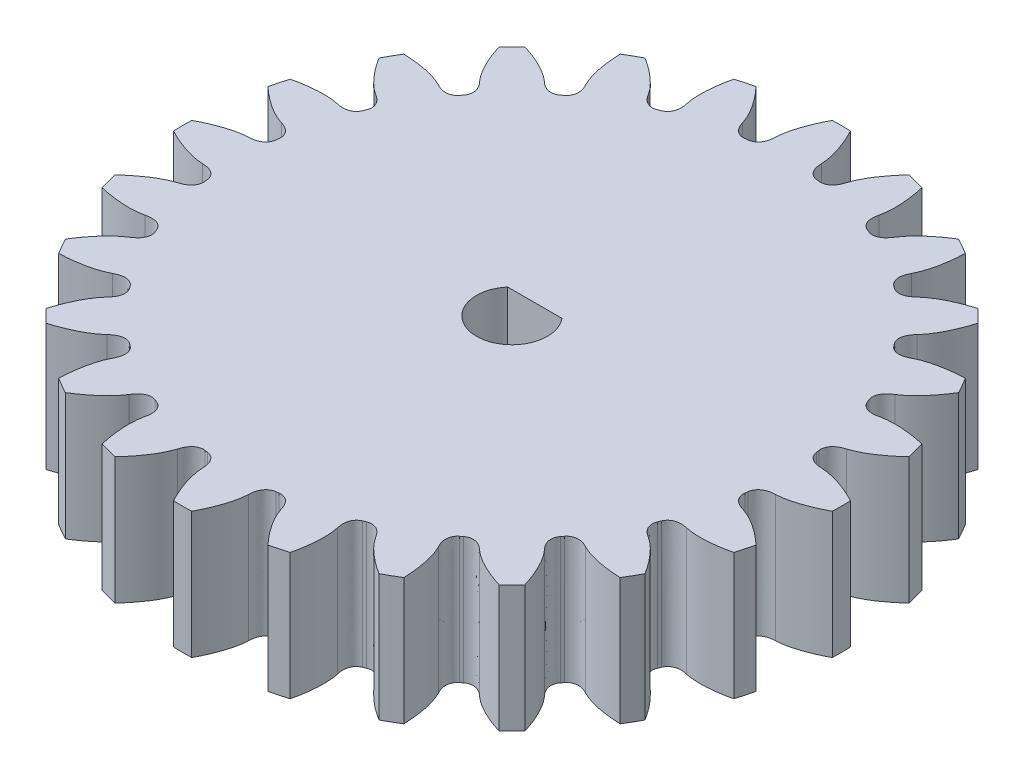
SolidWorks part; units mm, degrees
ref_plane "Спереди" through (0, 0, 0) normal (0, 0, 1) x (1, 0, 0)
ref_plane "Сверху" through (0, 0, 0) normal (0, 1, 0) x (1, 0, 0)
ref_plane "Справа" through (0, 0, 0) normal (1, 0, 0) x (0, 0, -1)
sketch "Эскиз1" plane through (0, 0, 0) normal (0, 1, 0) x (1, 0, 0)
  line L0 (-1.0724, 0.9) -> (1.0724, 0.9)
  arc A3 (-1.0724, 0.9) -> (1.0724, 0.9) centre (0, 0) ccw
  point P1 (0, -1.4)
  line B0 (-14.3, 0) -> (14.3, 0) construction
  line B1 (0, -14.3) -> (0, 14.3) construction
  arc B2 (0.3577, 12.9951) -> (-0.3577, 12.9951) centre (0, 0) ccw
  arc B3 (-1.346, 10.6654) -> (-1.4603, 10.6504) centre (0, 0) ccw
  arc B4 (-3.0178, 12.6449) -> (-3.7089, 12.4597) centre (0, 0) ccw
  arc B5 (-4.0605, 9.9536) -> (-4.1671, 9.9095) centre (0, 0) ccw
  arc B6 (-6.1877, 11.4329) -> (-6.8073, 11.0752) centre (0, 0) ccw
  arc B7 (-6.4984, 8.5635) -> (-6.5898, 8.4933) centre (0, 0) ccw
  arc B8 (-8.936, 9.4419) -> (-9.4419, 8.936) centre (0, 0) ccw
  arc B9 (-8.4933, 6.5898) -> (-8.5635, 6.4984) centre (0, 0) ccw
  arc B10 (-11.0752, 6.8073) -> (-11.4329, 6.1877) centre (0, 0) ccw
  arc B11 (-9.9095, 4.1671) -> (-9.9536, 4.0605) centre (0, 0) ccw
  arc B12 (-12.4597, 3.7089) -> (-12.6449, 3.0178) centre (0, 0) ccw
  arc B13 (-10.6504, 1.4603) -> (-10.6654, 1.346) centre (0, 0) ccw
  arc B14 (-12.9951, 0.3577) -> (-12.9951, -0.3577) centre (0, 0) ccw
  arc B15 (-10.6654, -1.346) -> (-10.6504, -1.4603) centre (0, 0) ccw
  arc B16 (-12.6449, -3.0178) -> (-12.4597, -3.7089) centre (0, 0) ccw
  arc B17 (-9.9536, -4.0605) -> (-9.9095, -4.1671) centre (0, 0) ccw
  arc B18 (-11.4329, -6.1877) -> (-11.0752, -6.8073) centre (0, 0) ccw
  arc B19 (-8.5635, -6.4984) -> (-8.4933, -6.5898) centre (0, 0) ccw
  arc B20 (-9.4419, -8.936) -> (-8.936, -9.4419) centre (0, 0) ccw
  arc B21 (-6.5898, -8.4933) -> (-6.4984, -8.5635) centre (0, 0) ccw
  arc B22 (-6.8073, -11.0752) -> (-6.1877, -11.4329) centre (0, 0) ccw
  arc B23 (-4.1671, -9.9095) -> (-4.0605, -9.9536) centre (0, 0) ccw
  arc B24 (-3.7089, -12.4597) -> (-3.0178, -12.6449) centre (0, 0) ccw
  arc B25 (-1.4603, -10.6504) -> (-1.346, -10.6654) centre (0, 0) ccw
  arc B26 (-0.3577, -12.9951) -> (0.3577, -12.9951) centre (0, 0) ccw
  arc B27 (1.346, -10.6654) -> (1.4603, -10.6504) centre (0, 0) ccw
  arc B28 (3.0178, -12.6449) -> (3.7089, -12.4597) centre (0, 0) ccw
  arc B29 (4.0605, -9.9536) -> (4.1671, -9.9095) centre (0, 0) ccw
  arc B30 (6.1877, -11.4329) -> (6.8073, -11.0752) centre (0, 0) ccw
  arc B31 (6.4984, -8.5635) -> (6.5898, -8.4933) centre (0, 0) ccw
  arc B32 (8.936, -9.4419) -> (9.4419, -8.936) centre (0, 0) ccw
  arc B33 (8.4933, -6.5898) -> (8.5635, -6.4984) centre (0, 0) ccw
  arc B34 (11.0752, -6.8073) -> (11.4329, -6.1877) centre (0, 0) ccw
  arc B35 (9.9095, -4.1671) -> (9.9536, -4.0605) centre (0, 0) ccw
  arc B36 (12.4597, -3.7089) -> (12.6449, -3.0178) centre (0, 0) ccw
  arc B37 (10.6504, -1.4603) -> (10.6654, -1.346) centre (0, 0) ccw
  arc B38 (12.9951, -0.3577) -> (12.9951, 0.3577) centre (0, 0) ccw
  arc B39 (10.6654, 1.346) -> (10.6504, 1.4603) centre (0, 0) ccw
  arc B40 (12.6449, 3.0178) -> (12.4597, 3.7089) centre (0, 0) ccw
  arc B41 (9.9536, 4.0605) -> (9.9095, 4.1671) centre (0, 0) ccw
  arc B42 (11.4329, 6.1877) -> (11.0752, 6.8073) centre (0, 0) ccw
  arc B43 (8.5635, 6.4984) -> (8.4933, 6.5898) centre (0, 0) ccw
  arc B44 (9.4419, 8.936) -> (8.936, 9.4419) centre (0, 0) ccw
  arc B45 (6.5898, 8.4933) -> (6.4984, 8.5635) centre (0, 0) ccw
  arc B46 (6.8073, 11.0752) -> (6.1877, 11.4329) centre (0, 0) ccw
  arc B47 (4.1671, 9.9095) -> (4.0605, 9.9536) centre (0, 0) ccw
  arc B48 (3.7089, 12.4597) -> (3.0178, 12.6449) centre (0, 0) ccw
  arc B49 (1.4603, 10.6504) -> (1.346, 10.6654) centre (0, 0) ccw
  circle B50 centre (0, 0) radius 12 construction
  spline B51 degree 3 poles (0.9058, 11.3017) (0.9058, 11.2304) (0.9138, 11.1608) (0.9299, 11.0929) (0.9396, 11.0522) (0.9513, 11.0113) (0.9676, 10.9727) (0.9799, 10.9437) (0.994, 10.915) (1.0107, 10.8883) (1.0248, 10.8656) (1.0406, 10.8436) (1.058, 10.8234) (1.0738, 10.805) (1.091, 10.7875) (1.1093, 10.7717) (1.1266, 10.7569) (1.1451, 10.7431) (1.1643, 10.7309) (1.1829, 10.7192) (1.2025, 10.7087) (1.2225, 10.6998) (1.2421, 10.6911) (1.2626, 10.6838) (1.2833, 10.678) (1.3038, 10.6723) (1.3247, 10.6681) (1.346, 10.6654) knots 0 0 0 0 1 1 1 2 2 2 3 3 3 4 4 4 5 5 5 6 6 6 7 7 7 8 8 8 9 9 9 9
  spline B52 degree 3 poles (-0.9058, 11.3017) (-0.9058, 11.2304) (-0.9138, 11.1608) (-0.9299, 11.0929) (-0.9396, 11.0522) (-0.9513, 11.0113) (-0.9676, 10.9727) (-0.9799, 10.9437) (-0.994, 10.915) (-1.0107, 10.8883) (-1.0248, 10.8656) (-1.0406, 10.8436) (-1.058, 10.8234) (-1.0738, 10.805) (-1.091, 10.7875) (-1.1093, 10.7717) (-1.1266, 10.7569) (-1.1451, 10.7431) (-1.1643, 10.7309) (-1.1829, 10.7192) (-1.2025, 10.7087) (-1.2225, 10.6998) (-1.2421, 10.6911) (-1.2626, 10.6838) (-1.2833, 10.678) (-1.3038, 10.6723) (-1.3247, 10.6681) (-1.346, 10.6654) knots 0 0 0 0 1 1 1 2 2 2 3 3 3 4 4 4 5 5 5 6 6 6 7 7 7 8 8 8 9 9 9 9
  spline B53 degree 3 poles (0.9058, 11.3017) (0.9032, 11.3642) (0.898, 11.4263) (0.8903, 11.4882) (0.8824, 11.551) (0.8712, 11.6136) (0.8589, 11.6757) (0.8463, 11.7389) (0.8314, 11.8016) (0.8153, 11.864) (0.7989, 11.9273) (0.7806, 11.9902) (0.7612, 12.0526) (0.7414, 12.116) (0.72, 12.179) (0.6975, 12.2415) (0.6746, 12.3049) (0.6503, 12.3678) (0.6249, 12.4303) (0.5991, 12.4937) (0.572, 12.5566) (0.5439, 12.6189) (0.5153, 12.6822) (0.4855, 12.745) (0.4547, 12.8073) (0.4235, 12.8704) (0.3912, 12.933) (0.3577, 12.9951) knots 0 0 0 0 1 1 1 2 2 2 3 3 3 4 4 4 5 5 5 6 6 6 7 7 7 8 8 8 9 9 9 9
  spline B54 degree 3 poles (-0.9058, 11.3017) (-0.9032, 11.3642) (-0.898, 11.4263) (-0.8903, 11.4882) (-0.8824, 11.551) (-0.8712, 11.6136) (-0.8589, 11.6757) (-0.8463, 11.7389) (-0.8314, 11.8016) (-0.8153, 11.864) (-0.7989, 11.9273) (-0.7806, 11.9902) (-0.7612, 12.0526) (-0.7414, 12.116) (-0.72, 12.179) (-0.6975, 12.2415) (-0.6746, 12.3049) (-0.6503, 12.3678) (-0.6249, 12.4303) (-0.5991, 12.4937) (-0.572, 12.5566) (-0.5439, 12.6189) (-0.5153, 12.6822) (-0.4855, 12.745) (-0.4547, 12.8073) (-0.4235, 12.8704) (-0.3912, 12.933) (-0.3577, 12.9951) knots 0 0 0 0 1 1 1 2 2 2 3 3 3 4 4 4 5 5 5 6 6 6 7 7 7 8 8 8 9 9 9 9
  spline B55 degree 3 poles (-2.0502, 11.151) (-2.0317, 11.0822) (-2.0059, 11.017) (-1.9728, 10.9556) (-1.9529, 10.9188) (-1.931, 10.8823) (-1.9053, 10.8493) (-1.886, 10.8244) (-1.8649, 10.8004) (-1.8419, 10.7789) (-1.8224, 10.7606) (-1.8014, 10.7435) (-1.7793, 10.7284) (-1.7594, 10.7148) (-1.7382, 10.7023) (-1.7164, 10.6918) (-1.6959, 10.6819) (-1.6745, 10.6734) (-1.6527, 10.6666) (-1.6318, 10.6601) (-1.6101, 10.655) (-1.5885, 10.6516) (-1.5672, 10.6483) (-1.5456, 10.6465) (-1.5241, 10.6463) (-1.5028, 10.6461) (-1.4816, 10.6475) (-1.4603, 10.6504) knots 0 0 0 0 1 1 1 2 2 2 3 3 3 4 4 4 5 5 5 6 6 6 7 7 7 8 8 8 9 9 9 9
  spline B56 degree 3 poles (-3.8, 10.6822) (-3.7815, 10.6133) (-3.7713, 10.544) (-3.7693, 10.4743) (-3.7681, 10.4325) (-3.7688, 10.3898) (-3.7746, 10.3484) (-3.7789, 10.3172) (-3.7852, 10.2858) (-3.7943, 10.2557) (-3.8021, 10.2302) (-3.8117, 10.2048) (-3.8232, 10.1807) (-3.8337, 10.1589) (-3.8458, 10.1376) (-3.8595, 10.1176) (-3.8723, 10.0988) (-3.8866, 10.0806) (-3.902, 10.0639) (-3.9169, 10.0478) (-3.9331, 10.0326) (-3.9502, 10.0188) (-3.9669, 10.0053) (-3.9848, 9.9929) (-4.0032, 9.982) (-4.0216, 9.9712) (-4.0406, 9.9618) (-4.0605, 9.9536) knots 0 0 0 0 1 1 1 2 2 2 3 3 3 4 4 4 5 5 5 6 6 6 7 7 7 8 8 8 9 9 9 9
  spline B57 degree 3 poles (-2.0502, 11.151) (-2.0689, 11.2107) (-2.09, 11.2694) (-2.1134, 11.3271) (-2.1373, 11.3858) (-2.1643, 11.4434) (-2.1923, 11.5002) (-2.2208, 11.5579) (-2.2514, 11.6147) (-2.2831, 11.6707) (-2.3153, 11.7276) (-2.3493, 11.7837) (-2.3842, 11.8389) (-2.4197, 11.8951) (-2.4567, 11.9503) (-2.4946, 12.0049) (-2.5331, 12.0602) (-2.5729, 12.1147) (-2.6136, 12.1685) (-2.6549, 12.223) (-2.6974, 12.2768) (-2.7407, 12.3297) (-2.7847, 12.3835) (-2.8297, 12.4364) (-2.8755, 12.4885) (-2.9221, 12.5415) (-2.9695, 12.5936) (-3.0178, 12.6449) knots 0 0 0 0 1 1 1 2 2 2 3 3 3 4 4 4 5 5 5 6 6 6 7 7 7 8 8 8 9 9 9 9
  spline B58 degree 3 poles (-3.8, 10.6822) (-3.8136, 10.7432) (-3.8247, 10.8046) (-3.8333, 10.8663) (-3.842, 10.929) (-3.8474, 10.9924) (-3.8515, 11.0556) (-3.8557, 11.1198) (-3.8576, 11.1843) (-3.8581, 11.2487) (-3.8587, 11.3141) (-3.8573, 11.3796) (-3.8547, 11.4449) (-3.852, 11.5113) (-3.8476, 11.5776) (-3.8421, 11.6438) (-3.8364, 11.711) (-3.8292, 11.7781) (-3.8208, 11.845) (-3.8123, 11.9129) (-3.8024, 11.9807) (-3.7914, 12.0482) (-3.7802, 12.1167) (-3.7676, 12.1851) (-3.754, 12.2532) (-3.7402, 12.3223) (-3.7251, 12.3911) (-3.7089, 12.4597) knots 0 0 0 0 1 1 1 2 2 2 3 3 3 4 4 4 5 5 5 6 6 6 7 7 7 8 8 8 9 9 9 9
  spline B59 degree 3 poles (-4.8664, 10.2404) (-4.8308, 10.1787) (-4.789, 10.1225) (-4.7411, 10.0717) (-4.7124, 10.0413) (-4.6817, 10.0117) (-4.6484, 9.9865) (-4.6233, 9.9675) (-4.5967, 9.9497) (-4.5689, 9.9349) (-4.5453, 9.9223) (-4.5206, 9.9111) (-4.4954, 9.9023) (-4.4726, 9.8943) (-4.4489, 9.8878) (-4.4252, 9.8833) (-4.4028, 9.879) (-4.3799, 9.8763) (-4.3571, 9.8754) (-4.3352, 9.8745) (-4.313, 9.8752) (-4.2912, 9.8776) (-4.2698, 9.8798) (-4.2484, 9.8837) (-4.2276, 9.8891) (-4.2071, 9.8944) (-4.1869, 9.9012) (-4.1671, 9.9095) knots 0 0 0 0 1 1 1 2 2 2 3 3 3 4 4 4 5 5 5 6 6 6 7 7 7 8 8 8 9 9 9 9
  spline B60 degree 3 poles (-6.4353, 9.3347) (-6.3996, 9.2729) (-6.3718, 9.2086) (-6.3518, 9.1418) (-6.3398, 9.1017) (-6.3295, 9.0604) (-6.3243, 9.0188) (-6.3204, 8.9876) (-6.3184, 8.9557) (-6.3194, 8.9242) (-6.3203, 8.8975) (-6.323, 8.8706) (-6.3279, 8.8443) (-6.3324, 8.8205) (-6.3386, 8.7968) (-6.3466, 8.7739) (-6.3541, 8.7524) (-6.3632, 8.7312) (-6.3738, 8.7111) (-6.384, 8.6917) (-6.3957, 8.6728) (-6.4086, 8.655) (-6.4213, 8.6377) (-6.4353, 8.6211) (-6.4504, 8.6058) (-6.4653, 8.5906) (-6.4813, 8.5765) (-6.4984, 8.5635) knots 0 0 0 0 1 1 1 2 2 2 3 3 3 4 4 4 5 5 5 6 6 6 7 7 7 8 8 8 9 9 9 9
  spline B61 degree 3 poles (-4.8664, 10.2404) (-4.8999, 10.2932) (-4.9355, 10.3445) (-4.9731, 10.3942) (-5.0113, 10.4447) (-5.0523, 10.4933) (-5.0941, 10.5409) (-5.1365, 10.5893) (-5.1808, 10.6362) (-5.2259, 10.6822) (-5.2718, 10.7288) (-5.319, 10.7741) (-5.3671, 10.8185) (-5.4159, 10.8635) (-5.4659, 10.9073) (-5.5167, 10.9502) (-5.5682, 10.9937) (-5.6207, 11.036) (-5.674, 11.0774) (-5.728, 11.1194) (-5.7829, 11.1603) (-5.8385, 11.2003) (-5.8949, 11.2408) (-5.9521, 11.2803) (-6.0098, 11.3188) (-6.0685, 11.3578) (-6.1278, 11.3959) (-6.1877, 11.4329) knots 0 0 0 0 1 1 1 2 2 2 3 3 3 4 4 4 5 5 5 6 6 6 7 7 7 8 8 8 9 9 9 9
  spline B62 degree 3 poles (-6.4353, 9.3347) (-6.4642, 9.3901) (-6.4908, 9.4465) (-6.5151, 9.5039) (-6.5397, 9.5623) (-6.5613, 9.622) (-6.5817, 9.6821) (-6.6024, 9.743) (-6.6209, 9.8048) (-6.638, 9.8669) (-6.6555, 9.9299) (-6.6711, 9.9935) (-6.6855, 10.0573) (-6.7001, 10.1221) (-6.713, 10.1873) (-6.7248, 10.2527) (-6.7367, 10.319) (-6.7471, 10.3857) (-6.7563, 10.4525) (-6.7657, 10.5203) (-6.7737, 10.5883) (-6.7805, 10.6564) (-6.7874, 10.7255) (-6.793, 10.7948) (-6.7974, 10.8641) (-6.8019, 10.9344) (-6.8053, 11.0047) (-6.8073, 11.0752) knots 0 0 0 0 1 1 1 2 2 2 3 3 3 4 4 4 5 5 5 6 6 6 7 7 7 8 8 8 9 9 9 9
  spline B63 degree 3 poles (-7.351, 8.632) (-7.3006, 8.5816) (-7.2457, 8.5381) (-7.1863, 8.5015) (-7.1507, 8.4795) (-7.1134, 8.4588) (-7.0747, 8.4431) (-7.0455, 8.4312) (-7.0152, 8.421) (-6.9845, 8.4138) (-6.9585, 8.4078) (-6.9318, 8.4034) (-6.9052, 8.4014) (-6.881, 8.3996) (-6.8565, 8.3994) (-6.8324, 8.4012) (-6.8097, 8.4029) (-6.7868, 8.4062) (-6.7646, 8.4112) (-6.7432, 8.416) (-6.7219, 8.4224) (-6.7015, 8.4304) (-6.6814, 8.4381) (-6.6618, 8.4474) (-6.6431, 8.4579) (-6.6246, 8.4684) (-6.6068, 8.4802) (-6.5898, 8.4933) knots 0 0 0 0 1 1 1 2 2 2 3 3 3 4 4 4 5 5 5 6 6 6 7 7 7 8 8 8 9 9 9 9
  spline B64 degree 3 poles (-8.632, 7.351) (-8.5816, 7.3006) (-8.5381, 7.2457) (-8.5015, 7.1863) (-8.4795, 7.1507) (-8.4588, 7.1134) (-8.4431, 7.0747) (-8.4312, 7.0455) (-8.421, 7.0152) (-8.4138, 6.9845) (-8.4078, 6.9585) (-8.4034, 6.9318) (-8.4014, 6.9052) (-8.3996, 6.881) (-8.3994, 6.8565) (-8.4012, 6.8324) (-8.4029, 6.8097) (-8.4062, 6.7868) (-8.4112, 6.7646) (-8.416, 6.7432) (-8.4224, 6.7219) (-8.4304, 6.7015) (-8.4381, 6.6814) (-8.4474, 6.6618) (-8.4579, 6.6431) (-8.4684, 6.6246) (-8.4802, 6.6068) (-8.4933, 6.5898) knots 0 0 0 0 1 1 1 2 2 2 3 3 3 4 4 4 5 5 5 6 6 6 7 7 7 8 8 8 9 9 9 9
  spline B65 degree 3 poles (-7.351, 8.632) (-7.3971, 8.6743) (-7.4447, 8.7146) (-7.4938, 8.7529) (-7.5438, 8.7918) (-7.596, 8.8281) (-7.6487, 8.8633) (-7.7022, 8.8991) (-7.7571, 8.9329) (-7.8126, 8.9656) (-7.869, 8.9988) (-7.9263, 9.0303) (-7.9843, 9.0607) (-8.0431, 9.0916) (-8.1027, 9.121) (-8.1628, 9.1492) (-8.2238, 9.1779) (-8.2855, 9.2052) (-8.3477, 9.2314) (-8.4107, 9.258) (-8.4744, 9.2833) (-8.5384, 9.3075) (-8.6033, 9.3321) (-8.6688, 9.3554) (-8.7346, 9.3776) (-8.8013, 9.4002) (-8.8684, 9.4216) (-8.936, 9.4419) knots 0 0 0 0 1 1 1 2 2 2 3 3 3 4 4 4 5 5 5 6 6 6 7 7 7 8 8 8 9 9 9 9
  spline B66 degree 3 poles (-8.632, 7.351) (-8.6743, 7.3971) (-8.7146, 7.4447) (-8.7529, 7.4938) (-8.7918, 7.5438) (-8.8281, 7.596) (-8.8633, 7.6487) (-8.8991, 7.7022) (-8.9329, 7.7571) (-8.9656, 7.8126) (-8.9988, 7.869) (-9.0303, 7.9263) (-9.0607, 7.9843) (-9.0916, 8.0431) (-9.121, 8.1027) (-9.1492, 8.1628) (-9.1779, 8.2238) (-9.2052, 8.2855) (-9.2314, 8.3477) (-9.258, 8.4107) (-9.2833, 8.4744) (-9.3075, 8.5384) (-9.3321, 8.6033) (-9.3554, 8.6688) (-9.3776, 8.7346) (-9.4002, 8.8013) (-9.4216, 8.8684) (-9.4419, 8.936) knots 0 0 0 0 1 1 1 2 2 2 3 3 3 4 4 4 5 5 5 6 6 6 7 7 7 8 8 8 9 9 9 9
  spline B67 degree 3 poles (-9.3347, 6.4353) (-9.2729, 6.3996) (-9.2086, 6.3718) (-9.1418, 6.3518) (-9.1017, 6.3398) (-9.0604, 6.3295) (-9.0188, 6.3243) (-8.9876, 6.3204) (-8.9557, 6.3184) (-8.9242, 6.3194) (-8.8975, 6.3203) (-8.8706, 6.323) (-8.8443, 6.3279) (-8.8205, 6.3324) (-8.7968, 6.3386) (-8.7739, 6.3466) (-8.7524, 6.3541) (-8.7312, 6.3632) (-8.7111, 6.3738) (-8.6917, 6.384) (-8.6728, 6.3957) (-8.655, 6.4086) (-8.6377, 6.4213) (-8.6211, 6.4353) (-8.6058, 6.4504) (-8.5906, 6.4653) (-8.5765, 6.4813) (-8.5635, 6.4984) knots 0 0 0 0 1 1 1 2 2 2 3 3 3 4 4 4 5 5 5 6 6 6 7 7 7 8 8 8 9 9 9 9
  spline B68 degree 3 poles (-10.2404, 4.8664) (-10.1787, 4.8308) (-10.1225, 4.789) (-10.0717, 4.7411) (-10.0413, 4.7124) (-10.0117, 4.6817) (-9.9865, 4.6484) (-9.9675, 4.6233) (-9.9497, 4.5967) (-9.9349, 4.5689) (-9.9223, 4.5453) (-9.9111, 4.5206) (-9.9023, 4.4954) (-9.8943, 4.4726) (-9.8878, 4.4489) (-9.8833, 4.4252) (-9.879, 4.4028) (-9.8763, 4.3799) (-9.8754, 4.3571) (-9.8745, 4.3352) (-9.8752, 4.313) (-9.8776, 4.2912) (-9.8798, 4.2698) (-9.8837, 4.2484) (-9.8891, 4.2276) (-9.8944, 4.2071) (-9.9012, 4.1869) (-9.9095, 4.1671) knots 0 0 0 0 1 1 1 2 2 2 3 3 3 4 4 4 5 5 5 6 6 6 7 7 7 8 8 8 9 9 9 9
  spline B69 degree 3 poles (-9.3347, 6.4353) (-9.3901, 6.4642) (-9.4465, 6.4908) (-9.5039, 6.5151) (-9.5623, 6.5397) (-9.622, 6.5613) (-9.6821, 6.5817) (-9.743, 6.6024) (-9.8048, 6.6209) (-9.8669, 6.638) (-9.9299, 6.6555) (-9.9935, 6.6711) (-10.0573, 6.6855) (-10.1221, 6.7001) (-10.1873, 6.713) (-10.2527, 6.7248) (-10.319, 6.7367) (-10.3857, 6.7471) (-10.4525, 6.7563) (-10.5203, 6.7657) (-10.5883, 6.7737) (-10.6564, 6.7805) (-10.7255, 6.7874) (-10.7948, 6.793) (-10.8641, 6.7974) (-10.9344, 6.8019) (-11.0047, 6.8053) (-11.0752, 6.8073) knots 0 0 0 0 1 1 1 2 2 2 3 3 3 4 4 4 5 5 5 6 6 6 7 7 7 8 8 8 9 9 9 9
  spline B70 degree 3 poles (-10.2404, 4.8664) (-10.2932, 4.8999) (-10.3445, 4.9355) (-10.3942, 4.9731) (-10.4447, 5.0113) (-10.4933, 5.0523) (-10.5409, 5.0941) (-10.5893, 5.1365) (-10.6362, 5.1808) (-10.6822, 5.2259) (-10.7288, 5.2718) (-10.7741, 5.319) (-10.8185, 5.3671) (-10.8635, 5.4159) (-10.9073, 5.4659) (-10.9502, 5.5167) (-10.9937, 5.5682) (-11.036, 5.6207) (-11.0774, 5.674) (-11.1194, 5.728) (-11.1603, 5.7829) (-11.2003, 5.8385) (-11.2408, 5.8949) (-11.2803, 5.9521) (-11.3188, 6.0098) (-11.3578, 6.0685) (-11.3959, 6.1278) (-11.4329, 6.1877) knots 0 0 0 0 1 1 1 2 2 2 3 3 3 4 4 4 5 5 5 6 6 6 7 7 7 8 8 8 9 9 9 9
  spline B71 degree 3 poles (-10.6822, 3.8) (-10.6133, 3.7815) (-10.544, 3.7713) (-10.4743, 3.7693) (-10.4325, 3.7681) (-10.3898, 3.7688) (-10.3484, 3.7746) (-10.3172, 3.7789) (-10.2858, 3.7852) (-10.2557, 3.7943) (-10.2302, 3.8021) (-10.2048, 3.8117) (-10.1807, 3.8232) (-10.1589, 3.8337) (-10.1376, 3.8458) (-10.1176, 3.8595) (-10.0988, 3.8723) (-10.0806, 3.8866) (-10.0639, 3.902) (-10.0478, 3.9169) (-10.0326, 3.9331) (-10.0188, 3.9502) (-10.0053, 3.9669) (-9.9929, 3.9848) (-9.982, 4.0032) (-9.9712, 4.0216) (-9.9618, 4.0406) (-9.9536, 4.0605) knots 0 0 0 0 1 1 1 2 2 2 3 3 3 4 4 4 5 5 5 6 6 6 7 7 7 8 8 8 9 9 9 9
  spline B72 degree 3 poles (-11.151, 2.0502) (-11.0822, 2.0317) (-11.017, 2.0059) (-10.9556, 1.9728) (-10.9188, 1.9529) (-10.8823, 1.931) (-10.8493, 1.9053) (-10.8244, 1.886) (-10.8004, 1.8649) (-10.7789, 1.8419) (-10.7606, 1.8224) (-10.7435, 1.8014) (-10.7284, 1.7793) (-10.7148, 1.7594) (-10.7023, 1.7382) (-10.6918, 1.7164) (-10.6819, 1.6959) (-10.6734, 1.6745) (-10.6666, 1.6527) (-10.6601, 1.6318) (-10.655, 1.6101) (-10.6516, 1.5885) (-10.6483, 1.5672) (-10.6465, 1.5456) (-10.6463, 1.5241) (-10.6461, 1.5028) (-10.6475, 1.4816) (-10.6504, 1.4603) knots 0 0 0 0 1 1 1 2 2 2 3 3 3 4 4 4 5 5 5 6 6 6 7 7 7 8 8 8 9 9 9 9
  spline B73 degree 3 poles (-10.6822, 3.8) (-10.7432, 3.8136) (-10.8046, 3.8247) (-10.8663, 3.8333) (-10.929, 3.842) (-10.9924, 3.8474) (-11.0556, 3.8515) (-11.1198, 3.8557) (-11.1843, 3.8576) (-11.2487, 3.8581) (-11.3141, 3.8587) (-11.3796, 3.8573) (-11.4449, 3.8547) (-11.5113, 3.852) (-11.5776, 3.8476) (-11.6438, 3.8421) (-11.711, 3.8364) (-11.7781, 3.8292) (-11.845, 3.8208) (-11.9129, 3.8123) (-11.9807, 3.8024) (-12.0482, 3.7914) (-12.1167, 3.7802) (-12.1851, 3.7676) (-12.2532, 3.754) (-12.3223, 3.7402) (-12.3911, 3.7251) (-12.4597, 3.7089) knots 0 0 0 0 1 1 1 2 2 2 3 3 3 4 4 4 5 5 5 6 6 6 7 7 7 8 8 8 9 9 9 9
  spline B74 degree 3 poles (-11.151, 2.0502) (-11.2107, 2.0689) (-11.2694, 2.09) (-11.3271, 2.1134) (-11.3858, 2.1373) (-11.4434, 2.1643) (-11.5002, 2.1923) (-11.5579, 2.2208) (-11.6147, 2.2514) (-11.6707, 2.2831) (-11.7276, 2.3153) (-11.7837, 2.3493) (-11.8389, 2.3842) (-11.8951, 2.4197) (-11.9503, 2.4567) (-12.0049, 2.4946) (-12.0602, 2.5331) (-12.1147, 2.5729) (-12.1685, 2.6136) (-12.223, 2.6549) (-12.2768, 2.6974) (-12.3297, 2.7407) (-12.3835, 2.7847) (-12.4364, 2.8297) (-12.4885, 2.8755) (-12.5415, 2.9221) (-12.5936, 2.9695) (-12.6449, 3.0178) knots 0 0 0 0 1 1 1 2 2 2 3 3 3 4 4 4 5 5 5 6 6 6 7 7 7 8 8 8 9 9 9 9
  spline B75 degree 3 poles (-11.3017, 0.9058) (-11.2304, 0.9058) (-11.1608, 0.9138) (-11.0929, 0.9299) (-11.0522, 0.9396) (-11.0113, 0.9513) (-10.9727, 0.9676) (-10.9437, 0.9799) (-10.915, 0.994) (-10.8883, 1.0107) (-10.8656, 1.0248) (-10.8436, 1.0406) (-10.8234, 1.058) (-10.805, 1.0738) (-10.7875, 1.091) (-10.7717, 1.1093) (-10.7569, 1.1266) (-10.7431, 1.1451) (-10.7309, 1.1643) (-10.7192, 1.1829) (-10.7087, 1.2025) (-10.6998, 1.2225) (-10.6911, 1.2421) (-10.6838, 1.2626) (-10.678, 1.2833) (-10.6723, 1.3038) (-10.6681, 1.3247) (-10.6654, 1.346) knots 0 0 0 0 1 1 1 2 2 2 3 3 3 4 4 4 5 5 5 6 6 6 7 7 7 8 8 8 9 9 9 9
  spline B76 degree 3 poles (-11.3017, -0.9058) (-11.2304, -0.9058) (-11.1608, -0.9138) (-11.0929, -0.9299) (-11.0522, -0.9396) (-11.0113, -0.9513) (-10.9727, -0.9676) (-10.9437, -0.9799) (-10.915, -0.994) (-10.8883, -1.0107) (-10.8656, -1.0248) (-10.8436, -1.0406) (-10.8234, -1.058) (-10.805, -1.0738) (-10.7875, -1.091) (-10.7717, -1.1093) (-10.7569, -1.1266) (-10.7431, -1.1451) (-10.7309, -1.1643) (-10.7192, -1.1829) (-10.7087, -1.2025) (-10.6998, -1.2225) (-10.6911, -1.2421) (-10.6838, -1.2626) (-10.678, -1.2833) (-10.6723, -1.3038) (-10.6681, -1.3247) (-10.6654, -1.346) knots 0 0 0 0 1 1 1 2 2 2 3 3 3 4 4 4 5 5 5 6 6 6 7 7 7 8 8 8 9 9 9 9
  spline B77 degree 3 poles (-11.3017, 0.9058) (-11.3642, 0.9032) (-11.4263, 0.898) (-11.4882, 0.8903) (-11.551, 0.8824) (-11.6136, 0.8712) (-11.6757, 0.8589) (-11.7389, 0.8463) (-11.8016, 0.8314) (-11.864, 0.8153) (-11.9273, 0.7989) (-11.9902, 0.7806) (-12.0526, 0.7612) (-12.116, 0.7414) (-12.179, 0.72) (-12.2415, 0.6975) (-12.3049, 0.6746) (-12.3678, 0.6503) (-12.4303, 0.6249) (-12.4937, 0.5991) (-12.5566, 0.572) (-12.6189, 0.5439) (-12.6822, 0.5153) (-12.745, 0.4855) (-12.8073, 0.4547) (-12.8704, 0.4235) (-12.933, 0.3912) (-12.9951, 0.3577) knots 0 0 0 0 1 1 1 2 2 2 3 3 3 4 4 4 5 5 5 6 6 6 7 7 7 8 8 8 9 9 9 9
  spline B78 degree 3 poles (-11.3017, -0.9058) (-11.3642, -0.9032) (-11.4263, -0.898) (-11.4882, -0.8903) (-11.551, -0.8824) (-11.6136, -0.8712) (-11.6757, -0.8589) (-11.7389, -0.8463) (-11.8016, -0.8314) (-11.864, -0.8153) (-11.9273, -0.7989) (-11.9902, -0.7806) (-12.0526, -0.7612) (-12.116, -0.7414) (-12.179, -0.72) (-12.2415, -0.6975) (-12.3049, -0.6746) (-12.3678, -0.6503) (-12.4303, -0.6249) (-12.4937, -0.5991) (-12.5566, -0.572) (-12.6189, -0.5439) (-12.6822, -0.5153) (-12.745, -0.4855) (-12.8073, -0.4547) (-12.8704, -0.4235) (-12.933, -0.3912) (-12.9951, -0.3577) knots 0 0 0 0 1 1 1 2 2 2 3 3 3 4 4 4 5 5 5 6 6 6 7 7 7 8 8 8 9 9 9 9
  spline B79 degree 3 poles (-11.151, -2.0502) (-11.0822, -2.0317) (-11.017, -2.0059) (-10.9556, -1.9728) (-10.9188, -1.9529) (-10.8823, -1.931) (-10.8493, -1.9053) (-10.8244, -1.886) (-10.8004, -1.8649) (-10.7789, -1.8419) (-10.7606, -1.8224) (-10.7435, -1.8014) (-10.7284, -1.7793) (-10.7148, -1.7594) (-10.7023, -1.7382) (-10.6918, -1.7164) (-10.6819, -1.6959) (-10.6734, -1.6745) (-10.6666, -1.6527) (-10.6601, -1.6318) (-10.655, -1.6101) (-10.6516, -1.5885) (-10.6483, -1.5672) (-10.6465, -1.5456) (-10.6463, -1.5241) (-10.6461, -1.5028) (-10.6475, -1.4816) (-10.6504, -1.4603) knots 0 0 0 0 1 1 1 2 2 2 3 3 3 4 4 4 5 5 5 6 6 6 7 7 7 8 8 8 9 9 9 9
  spline B80 degree 3 poles (-10.6822, -3.8) (-10.6133, -3.7815) (-10.544, -3.7713) (-10.4743, -3.7693) (-10.4325, -3.7681) (-10.3898, -3.7688) (-10.3484, -3.7746) (-10.3172, -3.7789) (-10.2858, -3.7852) (-10.2557, -3.7943) (-10.2302, -3.8021) (-10.2048, -3.8117) (-10.1807, -3.8232) (-10.1589, -3.8337) (-10.1376, -3.8458) (-10.1176, -3.8595) (-10.0988, -3.8723) (-10.0806, -3.8866) (-10.0639, -3.902) (-10.0478, -3.9169) (-10.0326, -3.9331) (-10.0188, -3.9502) (-10.0053, -3.9669) (-9.9929, -3.9848) (-9.982, -4.0032) (-9.9712, -4.0216) (-9.9618, -4.0406) (-9.9536, -4.0605) knots 0 0 0 0 1 1 1 2 2 2 3 3 3 4 4 4 5 5 5 6 6 6 7 7 7 8 8 8 9 9 9 9
  spline B81 degree 3 poles (-11.151, -2.0502) (-11.2107, -2.0689) (-11.2694, -2.09) (-11.3271, -2.1134) (-11.3858, -2.1373) (-11.4434, -2.1643) (-11.5002, -2.1923) (-11.5579, -2.2208) (-11.6147, -2.2514) (-11.6707, -2.2831) (-11.7276, -2.3153) (-11.7837, -2.3493) (-11.8389, -2.3842) (-11.8951, -2.4197) (-11.9503, -2.4567) (-12.0049, -2.4946) (-12.0602, -2.5331) (-12.1147, -2.5729) (-12.1685, -2.6136) (-12.223, -2.6549) (-12.2768, -2.6974) (-12.3297, -2.7407) (-12.3835, -2.7847) (-12.4364, -2.8297) (-12.4885, -2.8755) (-12.5415, -2.9221) (-12.5936, -2.9695) (-12.6449, -3.0178) knots 0 0 0 0 1 1 1 2 2 2 3 3 3 4 4 4 5 5 5 6 6 6 7 7 7 8 8 8 9 9 9 9
  spline B82 degree 3 poles (-10.6822, -3.8) (-10.7432, -3.8136) (-10.8046, -3.8247) (-10.8663, -3.8333) (-10.929, -3.842) (-10.9924, -3.8474) (-11.0556, -3.8515) (-11.1198, -3.8557) (-11.1843, -3.8576) (-11.2487, -3.8581) (-11.3141, -3.8587) (-11.3796, -3.8573) (-11.4449, -3.8547) (-11.5113, -3.852) (-11.5776, -3.8476) (-11.6438, -3.8421) (-11.711, -3.8364) (-11.7781, -3.8292) (-11.845, -3.8208) (-11.9129, -3.8123) (-11.9807, -3.8024) (-12.0482, -3.7914) (-12.1167, -3.7802) (-12.1851, -3.7676) (-12.2532, -3.754) (-12.3223, -3.7402) (-12.3911, -3.7251) (-12.4597, -3.7089) knots 0 0 0 0 1 1 1 2 2 2 3 3 3 4 4 4 5 5 5 6 6 6 7 7 7 8 8 8 9 9 9 9
  spline B83 degree 3 poles (-10.2404, -4.8664) (-10.1787, -4.8308) (-10.1225, -4.789) (-10.0717, -4.7411) (-10.0413, -4.7124) (-10.0117, -4.6817) (-9.9865, -4.6484) (-9.9675, -4.6233) (-9.9497, -4.5967) (-9.9349, -4.5689) (-9.9223, -4.5453) (-9.9111, -4.5206) (-9.9023, -4.4954) (-9.8943, -4.4726) (-9.8878, -4.4489) (-9.8833, -4.4252) (-9.879, -4.4028) (-9.8763, -4.3799) (-9.8754, -4.3571) (-9.8745, -4.3352) (-9.8752, -4.313) (-9.8776, -4.2912) (-9.8798, -4.2698) (-9.8837, -4.2484) (-9.8891, -4.2276) (-9.8944, -4.2071) (-9.9012, -4.1869) (-9.9095, -4.1671) knots 0 0 0 0 1 1 1 2 2 2 3 3 3 4 4 4 5 5 5 6 6 6 7 7 7 8 8 8 9 9 9 9
  spline B84 degree 3 poles (-9.3347, -6.4353) (-9.2729, -6.3996) (-9.2086, -6.3718) (-9.1418, -6.3518) (-9.1017, -6.3398) (-9.0604, -6.3295) (-9.0188, -6.3243) (-8.9876, -6.3204) (-8.9557, -6.3184) (-8.9242, -6.3194) (-8.8975, -6.3203) (-8.8706, -6.323) (-8.8443, -6.3279) (-8.8205, -6.3324) (-8.7968, -6.3386) (-8.7739, -6.3466) (-8.7524, -6.3541) (-8.7312, -6.3632) (-8.7111, -6.3738) (-8.6917, -6.384) (-8.6728, -6.3957) (-8.655, -6.4086) (-8.6377, -6.4213) (-8.6211, -6.4353) (-8.6058, -6.4504) (-8.5906, -6.4653) (-8.5765, -6.4813) (-8.5635, -6.4984) knots 0 0 0 0 1 1 1 2 2 2 3 3 3 4 4 4 5 5 5 6 6 6 7 7 7 8 8 8 9 9 9 9
  spline B85 degree 3 poles (-10.2404, -4.8664) (-10.2932, -4.8999) (-10.3445, -4.9355) (-10.3942, -4.9731) (-10.4447, -5.0113) (-10.4933, -5.0523) (-10.5409, -5.0941) (-10.5893, -5.1365) (-10.6362, -5.1808) (-10.6822, -5.2259) (-10.7288, -5.2718) (-10.7741, -5.319) (-10.8185, -5.3671) (-10.8635, -5.4159) (-10.9073, -5.4659) (-10.9502, -5.5167) (-10.9937, -5.5682) (-11.036, -5.6207) (-11.0774, -5.674) (-11.1194, -5.728) (-11.1603, -5.7829) (-11.2003, -5.8385) (-11.2408, -5.8949) (-11.2803, -5.9521) (-11.3188, -6.0098) (-11.3578, -6.0685) (-11.3959, -6.1278) (-11.4329, -6.1877) knots 0 0 0 0 1 1 1 2 2 2 3 3 3 4 4 4 5 5 5 6 6 6 7 7 7 8 8 8 9 9 9 9
  spline B86 degree 3 poles (-9.3347, -6.4353) (-9.3901, -6.4642) (-9.4465, -6.4908) (-9.5039, -6.5151) (-9.5623, -6.5397) (-9.622, -6.5613) (-9.6821, -6.5817) (-9.743, -6.6024) (-9.8048, -6.6209) (-9.8669, -6.638) (-9.9299, -6.6555) (-9.9935, -6.6711) (-10.0573, -6.6855) (-10.1221, -6.7001) (-10.1873, -6.713) (-10.2527, -6.7248) (-10.319, -6.7367) (-10.3857, -6.7471) (-10.4525, -6.7563) (-10.5203, -6.7657) (-10.5883, -6.7737) (-10.6564, -6.7805) (-10.7255, -6.7874) (-10.7948, -6.793) (-10.8641, -6.7974) (-10.9344, -6.8019) (-11.0047, -6.8053) (-11.0752, -6.8073) knots 0 0 0 0 1 1 1 2 2 2 3 3 3 4 4 4 5 5 5 6 6 6 7 7 7 8 8 8 9 9 9 9
  spline B87 degree 3 poles (-8.632, -7.351) (-8.5816, -7.3006) (-8.5381, -7.2457) (-8.5015, -7.1863) (-8.4795, -7.1507) (-8.4588, -7.1134) (-8.4431, -7.0747) (-8.4312, -7.0455) (-8.421, -7.0152) (-8.4138, -6.9845) (-8.4078, -6.9585) (-8.4034, -6.9318) (-8.4014, -6.9052) (-8.3996, -6.881) (-8.3994, -6.8565) (-8.4012, -6.8324) (-8.4029, -6.8097) (-8.4062, -6.7868) (-8.4112, -6.7646) (-8.416, -6.7432) (-8.4224, -6.7219) (-8.4304, -6.7015) (-8.4381, -6.6814) (-8.4474, -6.6618) (-8.4579, -6.6431) (-8.4684, -6.6246) (-8.4802, -6.6068) (-8.4933, -6.5898) knots 0 0 0 0 1 1 1 2 2 2 3 3 3 4 4 4 5 5 5 6 6 6 7 7 7 8 8 8 9 9 9 9
  spline B88 degree 3 poles (-7.351, -8.632) (-7.3006, -8.5816) (-7.2457, -8.5381) (-7.1863, -8.5015) (-7.1507, -8.4795) (-7.1134, -8.4588) (-7.0747, -8.4431) (-7.0455, -8.4312) (-7.0152, -8.421) (-6.9845, -8.4138) (-6.9585, -8.4078) (-6.9318, -8.4034) (-6.9052, -8.4014) (-6.881, -8.3996) (-6.8565, -8.3994) (-6.8324, -8.4012) (-6.8097, -8.4029) (-6.7868, -8.4062) (-6.7646, -8.4112) (-6.7432, -8.416) (-6.7219, -8.4224) (-6.7015, -8.4304) (-6.6814, -8.4381) (-6.6618, -8.4474) (-6.6431, -8.4579) (-6.6246, -8.4684) (-6.6068, -8.4802) (-6.5898, -8.4933) knots 0 0 0 0 1 1 1 2 2 2 3 3 3 4 4 4 5 5 5 6 6 6 7 7 7 8 8 8 9 9 9 9
  spline B89 degree 3 poles (-8.632, -7.351) (-8.6743, -7.3971) (-8.7146, -7.4447) (-8.7529, -7.4938) (-8.7918, -7.5438) (-8.8281, -7.596) (-8.8633, -7.6487) (-8.8991, -7.7022) (-8.9329, -7.7571) (-8.9656, -7.8126) (-8.9988, -7.869) (-9.0303, -7.9263) (-9.0607, -7.9843) (-9.0916, -8.0431) (-9.121, -8.1027) (-9.1492, -8.1628) (-9.1779, -8.2238) (-9.2052, -8.2855) (-9.2314, -8.3477) (-9.258, -8.4107) (-9.2833, -8.4744) (-9.3075, -8.5384) (-9.3321, -8.6033) (-9.3554, -8.6688) (-9.3776, -8.7346) (-9.4002, -8.8013) (-9.4216, -8.8684) (-9.4419, -8.936) knots 0 0 0 0 1 1 1 2 2 2 3 3 3 4 4 4 5 5 5 6 6 6 7 7 7 8 8 8 9 9 9 9
  spline B90 degree 3 poles (-7.351, -8.632) (-7.3971, -8.6743) (-7.4447, -8.7146) (-7.4938, -8.7529) (-7.5438, -8.7918) (-7.596, -8.8281) (-7.6487, -8.8633) (-7.7022, -8.8991) (-7.7571, -8.9329) (-7.8126, -8.9656) (-7.869, -8.9988) (-7.9263, -9.0303) (-7.9843, -9.0607) (-8.0431, -9.0916) (-8.1027, -9.121) (-8.1628, -9.1492) (-8.2238, -9.1779) (-8.2855, -9.2052) (-8.3477, -9.2314) (-8.4107, -9.258) (-8.4744, -9.2833) (-8.5384, -9.3075) (-8.6033, -9.3321) (-8.6688, -9.3554) (-8.7346, -9.3776) (-8.8013, -9.4002) (-8.8684, -9.4216) (-8.936, -9.4419) knots 0 0 0 0 1 1 1 2 2 2 3 3 3 4 4 4 5 5 5 6 6 6 7 7 7 8 8 8 9 9 9 9
  spline B91 degree 3 poles (-6.4353, -9.3347) (-6.3996, -9.2729) (-6.3718, -9.2086) (-6.3518, -9.1418) (-6.3398, -9.1017) (-6.3295, -9.0604) (-6.3243, -9.0188) (-6.3204, -8.9876) (-6.3184, -8.9557) (-6.3194, -8.9242) (-6.3203, -8.8975) (-6.323, -8.8706) (-6.3279, -8.8443) (-6.3324, -8.8205) (-6.3386, -8.7968) (-6.3466, -8.7739) (-6.3541, -8.7524) (-6.3632, -8.7312) (-6.3738, -8.7111) (-6.384, -8.6917) (-6.3957, -8.6728) (-6.4086, -8.655) (-6.4213, -8.6377) (-6.4353, -8.6211) (-6.4504, -8.6058) (-6.4653, -8.5906) (-6.4813, -8.5765) (-6.4984, -8.5635) knots 0 0 0 0 1 1 1 2 2 2 3 3 3 4 4 4 5 5 5 6 6 6 7 7 7 8 8 8 9 9 9 9
  spline B92 degree 3 poles (-4.8664, -10.2404) (-4.8308, -10.1787) (-4.789, -10.1225) (-4.7411, -10.0717) (-4.7124, -10.0413) (-4.6817, -10.0117) (-4.6484, -9.9865) (-4.6233, -9.9675) (-4.5967, -9.9497) (-4.5689, -9.9349) (-4.5453, -9.9223) (-4.5206, -9.9111) (-4.4954, -9.9023) (-4.4726, -9.8943) (-4.4489, -9.8878) (-4.4252, -9.8833) (-4.4028, -9.879) (-4.3799, -9.8763) (-4.3571, -9.8754) (-4.3352, -9.8745) (-4.313, -9.8752) (-4.2912, -9.8776) (-4.2698, -9.8798) (-4.2484, -9.8837) (-4.2276, -9.8891) (-4.2071, -9.8944) (-4.1869, -9.9012) (-4.1671, -9.9095) knots 0 0 0 0 1 1 1 2 2 2 3 3 3 4 4 4 5 5 5 6 6 6 7 7 7 8 8 8 9 9 9 9
  spline B93 degree 3 poles (-6.4353, -9.3347) (-6.4642, -9.3901) (-6.4908, -9.4465) (-6.5151, -9.5039) (-6.5397, -9.5623) (-6.5613, -9.622) (-6.5817, -9.6821) (-6.6024, -9.743) (-6.6209, -9.8048) (-6.638, -9.8669) (-6.6555, -9.9299) (-6.6711, -9.9935) (-6.6855, -10.0573) (-6.7001, -10.1221) (-6.713, -10.1873) (-6.7248, -10.2527) (-6.7367, -10.319) (-6.7471, -10.3857) (-6.7563, -10.4525) (-6.7657, -10.5203) (-6.7737, -10.5883) (-6.7805, -10.6564) (-6.7874, -10.7255) (-6.793, -10.7948) (-6.7974, -10.8641) (-6.8019, -10.9344) (-6.8053, -11.0047) (-6.8073, -11.0752) knots 0 0 0 0 1 1 1 2 2 2 3 3 3 4 4 4 5 5 5 6 6 6 7 7 7 8 8 8 9 9 9 9
  spline B94 degree 3 poles (-4.8664, -10.2404) (-4.8999, -10.2932) (-4.9355, -10.3445) (-4.9731, -10.3942) (-5.0113, -10.4447) (-5.0523, -10.4933) (-5.0941, -10.5409) (-5.1365, -10.5893) (-5.1808, -10.6362) (-5.2259, -10.6822) (-5.2718, -10.7288) (-5.319, -10.7741) (-5.3671, -10.8185) (-5.4159, -10.8635) (-5.4659, -10.9073) (-5.5167, -10.9502) (-5.5682, -10.9937) (-5.6207, -11.036) (-5.674, -11.0774) (-5.728, -11.1194) (-5.7829, -11.1603) (-5.8385, -11.2003) (-5.8949, -11.2408) (-5.9521, -11.2803) (-6.0098, -11.3188) (-6.0685, -11.3578) (-6.1278, -11.3959) (-6.1877, -11.4329) knots 0 0 0 0 1 1 1 2 2 2 3 3 3 4 4 4 5 5 5 6 6 6 7 7 7 8 8 8 9 9 9 9
  spline B95 degree 3 poles (-3.8, -10.6822) (-3.7815, -10.6133) (-3.7713, -10.544) (-3.7693, -10.4743) (-3.7681, -10.4325) (-3.7688, -10.3898) (-3.7746, -10.3484) (-3.7789, -10.3172) (-3.7852, -10.2858) (-3.7943, -10.2557) (-3.8021, -10.2302) (-3.8117, -10.2048) (-3.8232, -10.1807) (-3.8337, -10.1589) (-3.8458, -10.1376) (-3.8595, -10.1176) (-3.8723, -10.0988) (-3.8866, -10.0806) (-3.902, -10.0639) (-3.9169, -10.0478) (-3.9331, -10.0326) (-3.9502, -10.0188) (-3.9669, -10.0053) (-3.9848, -9.9929) (-4.0032, -9.982) (-4.0216, -9.9712) (-4.0406, -9.9618) (-4.0605, -9.9536) knots 0 0 0 0 1 1 1 2 2 2 3 3 3 4 4 4 5 5 5 6 6 6 7 7 7 8 8 8 9 9 9 9
  spline B96 degree 3 poles (-2.0502, -11.151) (-2.0317, -11.0822) (-2.0059, -11.017) (-1.9728, -10.9556) (-1.9529, -10.9188) (-1.931, -10.8823) (-1.9053, -10.8493) (-1.886, -10.8244) (-1.8649, -10.8004) (-1.8419, -10.7789) (-1.8224, -10.7606) (-1.8014, -10.7435) (-1.7793, -10.7284) (-1.7594, -10.7148) (-1.7382, -10.7023) (-1.7164, -10.6918) (-1.6959, -10.6819) (-1.6745, -10.6734) (-1.6527, -10.6666) (-1.6318, -10.6601) (-1.6101, -10.655) (-1.5885, -10.6516) (-1.5672, -10.6483) (-1.5456, -10.6465) (-1.5241, -10.6463) (-1.5028, -10.6461) (-1.4816, -10.6475) (-1.4603, -10.6504) knots 0 0 0 0 1 1 1 2 2 2 3 3 3 4 4 4 5 5 5 6 6 6 7 7 7 8 8 8 9 9 9 9
  spline B97 degree 3 poles (-3.8, -10.6822) (-3.8136, -10.7432) (-3.8247, -10.8046) (-3.8333, -10.8663) (-3.842, -10.929) (-3.8474, -10.9924) (-3.8515, -11.0556) (-3.8557, -11.1198) (-3.8576, -11.1843) (-3.8581, -11.2487) (-3.8587, -11.3141) (-3.8573, -11.3796) (-3.8547, -11.4449) (-3.852, -11.5113) (-3.8476, -11.5776) (-3.8421, -11.6438) (-3.8364, -11.711) (-3.8292, -11.7781) (-3.8208, -11.845) (-3.8123, -11.9129) (-3.8024, -11.9807) (-3.7914, -12.0482) (-3.7802, -12.1167) (-3.7676, -12.1851) (-3.754, -12.2532) (-3.7402, -12.3223) (-3.7251, -12.3911) (-3.7089, -12.4597) knots 0 0 0 0 1 1 1 2 2 2 3 3 3 4 4 4 5 5 5 6 6 6 7 7 7 8 8 8 9 9 9 9
  spline B98 degree 3 poles (-2.0502, -11.151) (-2.0689, -11.2107) (-2.09, -11.2694) (-2.1134, -11.3271) (-2.1373, -11.3858) (-2.1643, -11.4434) (-2.1923, -11.5002) (-2.2208, -11.5579) (-2.2514, -11.6147) (-2.2831, -11.6707) (-2.3153, -11.7276) (-2.3493, -11.7837) (-2.3842, -11.8389) (-2.4197, -11.8951) (-2.4567, -11.9503) (-2.4946, -12.0049) (-2.5331, -12.0602) (-2.5729, -12.1147) (-2.6136, -12.1685) (-2.6549, -12.223) (-2.6974, -12.2768) (-2.7407, -12.3297) (-2.7847, -12.3835) (-2.8297, -12.4364) (-2.8755, -12.4885) (-2.9221, -12.5415) (-2.9695, -12.5936) (-3.0178, -12.6449) knots 0 0 0 0 1 1 1 2 2 2 3 3 3 4 4 4 5 5 5 6 6 6 7 7 7 8 8 8 9 9 9 9
  spline B99 degree 3 poles (-0.9058, -11.3017) (-0.9058, -11.2304) (-0.9138, -11.1608) (-0.9299, -11.0929) (-0.9396, -11.0522) (-0.9513, -11.0113) (-0.9676, -10.9727) (-0.9799, -10.9437) (-0.994, -10.915) (-1.0107, -10.8883) (-1.0248, -10.8656) (-1.0406, -10.8436) (-1.058, -10.8234) (-1.0738, -10.805) (-1.091, -10.7875) (-1.1093, -10.7717) (-1.1266, -10.7569) (-1.1451, -10.7431) (-1.1643, -10.7309) (-1.1829, -10.7192) (-1.2025, -10.7087) (-1.2225, -10.6998) (-1.2421, -10.6911) (-1.2626, -10.6838) (-1.2833, -10.678) (-1.3038, -10.6723) (-1.3247, -10.6681) (-1.346, -10.6654) knots 0 0 0 0 1 1 1 2 2 2 3 3 3 4 4 4 5 5 5 6 6 6 7 7 7 8 8 8 9 9 9 9
  spline B100 degree 3 poles (0.9058, -11.3017) (0.9058, -11.2304) (0.9138, -11.1608) (0.9299, -11.0929) (0.9396, -11.0522) (0.9513, -11.0113) (0.9676, -10.9727) (0.9799, -10.9437) (0.994, -10.915) (1.0107, -10.8883) (1.0248, -10.8656) (1.0406, -10.8436) (1.058, -10.8234) (1.0738, -10.805) (1.091, -10.7875) (1.1093, -10.7717) (1.1266, -10.7569) (1.1451, -10.7431) (1.1643, -10.7309) (1.1829, -10.7192) (1.2025, -10.7087) (1.2225, -10.6998) (1.2421, -10.6911) (1.2626, -10.6838) (1.2833, -10.678) (1.3038, -10.6723) (1.3247, -10.6681) (1.346, -10.6654) knots 0 0 0 0 1 1 1 2 2 2 3 3 3 4 4 4 5 5 5 6 6 6 7 7 7 8 8 8 9 9 9 9
  spline B101 degree 3 poles (-0.9058, -11.3017) (-0.9032, -11.3642) (-0.898, -11.4263) (-0.8903, -11.4882) (-0.8824, -11.551) (-0.8712, -11.6136) (-0.8589, -11.6757) (-0.8463, -11.7389) (-0.8314, -11.8016) (-0.8153, -11.864) (-0.7989, -11.9273) (-0.7806, -11.9902) (-0.7612, -12.0526) (-0.7414, -12.116) (-0.72, -12.179) (-0.6975, -12.2415) (-0.6746, -12.3049) (-0.6503, -12.3678) (-0.6249, -12.4303) (-0.5991, -12.4937) (-0.572, -12.5566) (-0.5439, -12.6189) (-0.5153, -12.6822) (-0.4855, -12.745) (-0.4547, -12.8073) (-0.4235, -12.8704) (-0.3912, -12.933) (-0.3577, -12.9951) knots 0 0 0 0 1 1 1 2 2 2 3 3 3 4 4 4 5 5 5 6 6 6 7 7 7 8 8 8 9 9 9 9
  spline B102 degree 3 poles (0.9058, -11.3017) (0.9032, -11.3642) (0.898, -11.4263) (0.8903, -11.4882) (0.8824, -11.551) (0.8712, -11.6136) (0.8589, -11.6757) (0.8463, -11.7389) (0.8314, -11.8016) (0.8153, -11.864) (0.7989, -11.9273) (0.7806, -11.9902) (0.7612, -12.0526) (0.7414, -12.116) (0.72, -12.179) (0.6975, -12.2415) (0.6746, -12.3049) (0.6503, -12.3678) (0.6249, -12.4303) (0.5991, -12.4937) (0.572, -12.5566) (0.5439, -12.6189) (0.5153, -12.6822) (0.4855, -12.745) (0.4547, -12.8073) (0.4235, -12.8704) (0.3912, -12.933) (0.3577, -12.9951) knots 0 0 0 0 1 1 1 2 2 2 3 3 3 4 4 4 5 5 5 6 6 6 7 7 7 8 8 8 9 9 9 9
  spline B103 degree 3 poles (2.0502, -11.151) (2.0317, -11.0822) (2.0059, -11.017) (1.9728, -10.9556) (1.9529, -10.9188) (1.931, -10.8823) (1.9053, -10.8493) (1.886, -10.8244) (1.8649, -10.8004) (1.8419, -10.7789) (1.8224, -10.7606) (1.8014, -10.7435) (1.7793, -10.7284) (1.7594, -10.7148) (1.7382, -10.7023) (1.7164, -10.6918) (1.6959, -10.6819) (1.6745, -10.6734) (1.6527, -10.6666) (1.6318, -10.6601) (1.6101, -10.655) (1.5885, -10.6516) (1.5672, -10.6483) (1.5456, -10.6465) (1.5241, -10.6463) (1.5028, -10.6461) (1.4816, -10.6475) (1.4603, -10.6504) knots 0 0 0 0 1 1 1 2 2 2 3 3 3 4 4 4 5 5 5 6 6 6 7 7 7 8 8 8 9 9 9 9
  spline B104 degree 3 poles (3.8, -10.6822) (3.7815, -10.6133) (3.7713, -10.544) (3.7693, -10.4743) (3.7681, -10.4325) (3.7688, -10.3898) (3.7746, -10.3484) (3.7789, -10.3172) (3.7852, -10.2858) (3.7943, -10.2557) (3.8021, -10.2302) (3.8117, -10.2048) (3.8232, -10.1807) (3.8337, -10.1589) (3.8458, -10.1376) (3.8595, -10.1176) (3.8723, -10.0988) (3.8866, -10.0806) (3.902, -10.0639) (3.9169, -10.0478) (3.9331, -10.0326) (3.9502, -10.0188) (3.9669, -10.0053) (3.9848, -9.9929) (4.0032, -9.982) (4.0216, -9.9712) (4.0406, -9.9618) (4.0605, -9.9536) knots 0 0 0 0 1 1 1 2 2 2 3 3 3 4 4 4 5 5 5 6 6 6 7 7 7 8 8 8 9 9 9 9
  spline B105 degree 3 poles (2.0502, -11.151) (2.0689, -11.2107) (2.09, -11.2694) (2.1134, -11.3271) (2.1373, -11.3858) (2.1643, -11.4434) (2.1923, -11.5002) (2.2208, -11.5579) (2.2514, -11.6147) (2.2831, -11.6707) (2.3153, -11.7276) (2.3493, -11.7837) (2.3842, -11.8389) (2.4197, -11.8951) (2.4567, -11.9503) (2.4946, -12.0049) (2.5331, -12.0602) (2.5729, -12.1147) (2.6136, -12.1685) (2.6549, -12.223) (2.6974, -12.2768) (2.7407, -12.3297) (2.7847, -12.3835) (2.8297, -12.4364) (2.8755, -12.4885) (2.9221, -12.5415) (2.9695, -12.5936) (3.0178, -12.6449) knots 0 0 0 0 1 1 1 2 2 2 3 3 3 4 4 4 5 5 5 6 6 6 7 7 7 8 8 8 9 9 9 9
  spline B106 degree 3 poles (3.8, -10.6822) (3.8136, -10.7432) (3.8247, -10.8046) (3.8333, -10.8663) (3.842, -10.929) (3.8474, -10.9924) (3.8515, -11.0556) (3.8557, -11.1198) (3.8576, -11.1843) (3.8581, -11.2487) (3.8587, -11.3141) (3.8573, -11.3796) (3.8547, -11.4449) (3.852, -11.5113) (3.8476, -11.5776) (3.8421, -11.6438) (3.8364, -11.711) (3.8292, -11.7781) (3.8208, -11.845) (3.8123, -11.9129) (3.8024, -11.9807) (3.7914, -12.0482) (3.7802, -12.1167) (3.7676, -12.1851) (3.754, -12.2532) (3.7402, -12.3223) (3.7251, -12.3911) (3.7089, -12.4597) knots 0 0 0 0 1 1 1 2 2 2 3 3 3 4 4 4 5 5 5 6 6 6 7 7 7 8 8 8 9 9 9 9
  spline B107 degree 3 poles (4.8664, -10.2404) (4.8308, -10.1787) (4.789, -10.1225) (4.7411, -10.0717) (4.7124, -10.0413) (4.6817, -10.0117) (4.6484, -9.9865) (4.6233, -9.9675) (4.5967, -9.9497) (4.5689, -9.9349) (4.5453, -9.9223) (4.5206, -9.9111) (4.4954, -9.9023) (4.4726, -9.8943) (4.4489, -9.8878) (4.4252, -9.8833) (4.4028, -9.879) (4.3799, -9.8763) (4.3571, -9.8754) (4.3352, -9.8745) (4.313, -9.8752) (4.2912, -9.8776) (4.2698, -9.8798) (4.2484, -9.8837) (4.2276, -9.8891) (4.2071, -9.8944) (4.1869, -9.9012) (4.1671, -9.9095) knots 0 0 0 0 1 1 1 2 2 2 3 3 3 4 4 4 5 5 5 6 6 6 7 7 7 8 8 8 9 9 9 9
  spline B108 degree 3 poles (6.4353, -9.3347) (6.3996, -9.2729) (6.3718, -9.2086) (6.3518, -9.1418) (6.3398, -9.1017) (6.3295, -9.0604) (6.3243, -9.0188) (6.3204, -8.9876) (6.3184, -8.9557) (6.3194, -8.9242) (6.3203, -8.8975) (6.323, -8.8706) (6.3279, -8.8443) (6.3324, -8.8205) (6.3386, -8.7968) (6.3466, -8.7739) (6.3541, -8.7524) (6.3632, -8.7312) (6.3738, -8.7111) (6.384, -8.6917) (6.3957, -8.6728) (6.4086, -8.655) (6.4213, -8.6377) (6.4353, -8.6211) (6.4504, -8.6058) (6.4653, -8.5906) (6.4813, -8.5765) (6.4984, -8.5635) knots 0 0 0 0 1 1 1 2 2 2 3 3 3 4 4 4 5 5 5 6 6 6 7 7 7 8 8 8 9 9 9 9
  spline B109 degree 3 poles (4.8664, -10.2404) (4.8999, -10.2932) (4.9355, -10.3445) (4.9731, -10.3942) (5.0113, -10.4447) (5.0523, -10.4933) (5.0941, -10.5409) (5.1365, -10.5893) (5.1808, -10.6362) (5.2259, -10.6822) (5.2718, -10.7288) (5.319, -10.7741) (5.3671, -10.8185) (5.4159, -10.8635) (5.4659, -10.9073) (5.5167, -10.9502) (5.5682, -10.9937) (5.6207, -11.036) (5.674, -11.0774) (5.728, -11.1194) (5.7829, -11.1603) (5.8385, -11.2003) (5.8949, -11.2408) (5.9521, -11.2803) (6.0098, -11.3188) (6.0685, -11.3578) (6.1278, -11.3959) (6.1877, -11.4329) knots 0 0 0 0 1 1 1 2 2 2 3 3 3 4 4 4 5 5 5 6 6 6 7 7 7 8 8 8 9 9 9 9
  spline B110 degree 3 poles (6.4353, -9.3347) (6.4642, -9.3901) (6.4908, -9.4465) (6.5151, -9.5039) (6.5397, -9.5623) (6.5613, -9.622) (6.5817, -9.6821) (6.6024, -9.743) (6.6209, -9.8048) (6.638, -9.8669) (6.6555, -9.9299) (6.6711, -9.9935) (6.6855, -10.0573) (6.7001, -10.1221) (6.713, -10.1873) (6.7248, -10.2527) (6.7367, -10.319) (6.7471, -10.3857) (6.7563, -10.4525) (6.7657, -10.5203) (6.7737, -10.5883) (6.7805, -10.6564) (6.7874, -10.7255) (6.793, -10.7948) (6.7974, -10.8641) (6.8019, -10.9344) (6.8053, -11.0047) (6.8073, -11.0752) knots 0 0 0 0 1 1 1 2 2 2 3 3 3 4 4 4 5 5 5 6 6 6 7 7 7 8 8 8 9 9 9 9
  spline B111 degree 3 poles (7.351, -8.632) (7.3006, -8.5816) (7.2457, -8.5381) (7.1863, -8.5015) (7.1507, -8.4795) (7.1134, -8.4588) (7.0747, -8.4431) (7.0455, -8.4312) (7.0152, -8.421) (6.9845, -8.4138) (6.9585, -8.4078) (6.9318, -8.4034) (6.9052, -8.4014) (6.881, -8.3996) (6.8565, -8.3994) (6.8324, -8.4012) (6.8097, -8.4029) (6.7868, -8.4062) (6.7646, -8.4112) (6.7432, -8.416) (6.7219, -8.4224) (6.7015, -8.4304) (6.6814, -8.4381) (6.6618, -8.4474) (6.6431, -8.4579) (6.6246, -8.4684) (6.6068, -8.4802) (6.5898, -8.4933) knots 0 0 0 0 1 1 1 2 2 2 3 3 3 4 4 4 5 5 5 6 6 6 7 7 7 8 8 8 9 9 9 9
  spline B112 degree 3 poles (8.632, -7.351) (8.5816, -7.3006) (8.5381, -7.2457) (8.5015, -7.1863) (8.4795, -7.1507) (8.4588, -7.1134) (8.4431, -7.0747) (8.4312, -7.0455) (8.421, -7.0152) (8.4138, -6.9845) (8.4078, -6.9585) (8.4034, -6.9318) (8.4014, -6.9052) (8.3996, -6.881) (8.3994, -6.8565) (8.4012, -6.8324) (8.4029, -6.8097) (8.4062, -6.7868) (8.4112, -6.7646) (8.416, -6.7432) (8.4224, -6.7219) (8.4304, -6.7015) (8.4381, -6.6814) (8.4474, -6.6618) (8.4579, -6.6431) (8.4684, -6.6246) (8.4802, -6.6068) (8.4933, -6.5898) knots 0 0 0 0 1 1 1 2 2 2 3 3 3 4 4 4 5 5 5 6 6 6 7 7 7 8 8 8 9 9 9 9
  spline B113 degree 3 poles (7.351, -8.632) (7.3971, -8.6743) (7.4447, -8.7146) (7.4938, -8.7529) (7.5438, -8.7918) (7.596, -8.8281) (7.6487, -8.8633) (7.7022, -8.8991) (7.7571, -8.9329) (7.8126, -8.9656) (7.869, -8.9988) (7.9263, -9.0303) (7.9843, -9.0607) (8.0431, -9.0916) (8.1027, -9.121) (8.1628, -9.1492) (8.2238, -9.1779) (8.2855, -9.2052) (8.3477, -9.2314) (8.4107, -9.258) (8.4744, -9.2833) (8.5384, -9.3075) (8.6033, -9.3321) (8.6688, -9.3554) (8.7346, -9.3776) (8.8013, -9.4002) (8.8684, -9.4216) (8.936, -9.4419) knots 0 0 0 0 1 1 1 2 2 2 3 3 3 4 4 4 5 5 5 6 6 6 7 7 7 8 8 8 9 9 9 9
  spline B114 degree 3 poles (8.632, -7.351) (8.6743, -7.3971) (8.7146, -7.4447) (8.7529, -7.4938) (8.7918, -7.5438) (8.8281, -7.596) (8.8633, -7.6487) (8.8991, -7.7022) (8.9329, -7.7571) (8.9656, -7.8126) (8.9988, -7.869) (9.0303, -7.9263) (9.0607, -7.9843) (9.0916, -8.0431) (9.121, -8.1027) (9.1492, -8.1628) (9.1779, -8.2238) (9.2052, -8.2855) (9.2314, -8.3477) (9.258, -8.4107) (9.2833, -8.4744) (9.3075, -8.5384) (9.3321, -8.6033) (9.3554, -8.6688) (9.3776, -8.7346) (9.4002, -8.8013) (9.4216, -8.8684) (9.4419, -8.936) knots 0 0 0 0 1 1 1 2 2 2 3 3 3 4 4 4 5 5 5 6 6 6 7 7 7 8 8 8 9 9 9 9
  spline B115 degree 3 poles (9.3347, -6.4353) (9.2729, -6.3996) (9.2086, -6.3718) (9.1418, -6.3518) (9.1017, -6.3398) (9.0604, -6.3295) (9.0188, -6.3243) (8.9876, -6.3204) (8.9557, -6.3184) (8.9242, -6.3194) (8.8975, -6.3203) (8.8706, -6.323) (8.8443, -6.3279) (8.8205, -6.3324) (8.7968, -6.3386) (8.7739, -6.3466) (8.7524, -6.3541) (8.7312, -6.3632) (8.7111, -6.3738) (8.6917, -6.384) (8.6728, -6.3957) (8.655, -6.4086) (8.6377, -6.4213) (8.6211, -6.4353) (8.6058, -6.4504) (8.5906, -6.4653) (8.5765, -6.4813) (8.5635, -6.4984) knots 0 0 0 0 1 1 1 2 2 2 3 3 3 4 4 4 5 5 5 6 6 6 7 7 7 8 8 8 9 9 9 9
  spline B116 degree 3 poles (10.2404, -4.8664) (10.1787, -4.8308) (10.1225, -4.789) (10.0717, -4.7411) (10.0413, -4.7124) (10.0117, -4.6817) (9.9865, -4.6484) (9.9675, -4.6233) (9.9497, -4.5967) (9.9349, -4.5689) (9.9223, -4.5453) (9.9111, -4.5206) (9.9023, -4.4954) (9.8943, -4.4726) (9.8878, -4.4489) (9.8833, -4.4252) (9.879, -4.4028) (9.8763, -4.3799) (9.8754, -4.3571) (9.8745, -4.3352) (9.8752, -4.313) (9.8776, -4.2912) (9.8798, -4.2698) (9.8837, -4.2484) (9.8891, -4.2276) (9.8944, -4.2071) (9.9012, -4.1869) (9.9095, -4.1671) knots 0 0 0 0 1 1 1 2 2 2 3 3 3 4 4 4 5 5 5 6 6 6 7 7 7 8 8 8 9 9 9 9
  spline B117 degree 3 poles (9.3347, -6.4353) (9.3901, -6.4642) (9.4465, -6.4908) (9.5039, -6.5151) (9.5623, -6.5397) (9.622, -6.5613) (9.6821, -6.5817) (9.743, -6.6024) (9.8048, -6.6209) (9.8669, -6.638) (9.9299, -6.6555) (9.9935, -6.6711) (10.0573, -6.6855) (10.1221, -6.7001) (10.1873, -6.713) (10.2527, -6.7248) (10.319, -6.7367) (10.3857, -6.7471) (10.4525, -6.7563) (10.5203, -6.7657) (10.5883, -6.7737) (10.6564, -6.7805) (10.7255, -6.7874) (10.7948, -6.793) (10.8641, -6.7974) (10.9344, -6.8019) (11.0047, -6.8053) (11.0752, -6.8073) knots 0 0 0 0 1 1 1 2 2 2 3 3 3 4 4 4 5 5 5 6 6 6 7 7 7 8 8 8 9 9 9 9
  spline B118 degree 3 poles (10.2404, -4.8664) (10.2932, -4.8999) (10.3445, -4.9355) (10.3942, -4.9731) (10.4447, -5.0113) (10.4933, -5.0523) (10.5409, -5.0941) (10.5893, -5.1365) (10.6362, -5.1808) (10.6822, -5.2259) (10.7288, -5.2718) (10.7741, -5.319) (10.8185, -5.3671) (10.8635, -5.4159) (10.9073, -5.4659) (10.9502, -5.5167) (10.9937, -5.5682) (11.036, -5.6207) (11.0774, -5.674) (11.1194, -5.728) (11.1603, -5.7829) (11.2003, -5.8385) (11.2408, -5.8949) (11.2803, -5.9521) (11.3188, -6.0098) (11.3578, -6.0685) (11.3959, -6.1278) (11.4329, -6.1877) knots 0 0 0 0 1 1 1 2 2 2 3 3 3 4 4 4 5 5 5 6 6 6 7 7 7 8 8 8 9 9 9 9
  spline B119 degree 3 poles (10.6822, -3.8) (10.6133, -3.7815) (10.544, -3.7713) (10.4743, -3.7693) (10.4325, -3.7681) (10.3898, -3.7688) (10.3484, -3.7746) (10.3172, -3.7789) (10.2858, -3.7852) (10.2557, -3.7943) (10.2302, -3.8021) (10.2048, -3.8117) (10.1807, -3.8232) (10.1589, -3.8337) (10.1376, -3.8458) (10.1176, -3.8595) (10.0988, -3.8723) (10.0806, -3.8866) (10.0639, -3.902) (10.0478, -3.9169) (10.0326, -3.9331) (10.0188, -3.9502) (10.0053, -3.9669) (9.9929, -3.9848) (9.982, -4.0032) (9.9712, -4.0216) (9.9618, -4.0406) (9.9536, -4.0605) knots 0 0 0 0 1 1 1 2 2 2 3 3 3 4 4 4 5 5 5 6 6 6 7 7 7 8 8 8 9 9 9 9
  spline B120 degree 3 poles (11.151, -2.0502) (11.0822, -2.0317) (11.017, -2.0059) (10.9556, -1.9728) (10.9188, -1.9529) (10.8823, -1.931) (10.8493, -1.9053) (10.8244, -1.886) (10.8004, -1.8649) (10.7789, -1.8419) (10.7606, -1.8224) (10.7435, -1.8014) (10.7284, -1.7793) (10.7148, -1.7594) (10.7023, -1.7382) (10.6918, -1.7164) (10.6819, -1.6959) (10.6734, -1.6745) (10.6666, -1.6527) (10.6601, -1.6318) (10.655, -1.6101) (10.6516, -1.5885) (10.6483, -1.5672) (10.6465, -1.5456) (10.6463, -1.5241) (10.6461, -1.5028) (10.6475, -1.4816) (10.6504, -1.4603) knots 0 0 0 0 1 1 1 2 2 2 3 3 3 4 4 4 5 5 5 6 6 6 7 7 7 8 8 8 9 9 9 9
  spline B121 degree 3 poles (10.6822, -3.8) (10.7432, -3.8136) (10.8046, -3.8247) (10.8663, -3.8333) (10.929, -3.842) (10.9924, -3.8474) (11.0556, -3.8515) (11.1198, -3.8557) (11.1843, -3.8576) (11.2487, -3.8581) (11.3141, -3.8587) (11.3796, -3.8573) (11.4449, -3.8547) (11.5113, -3.852) (11.5776, -3.8476) (11.6438, -3.8421) (11.711, -3.8364) (11.7781, -3.8292) (11.845, -3.8208) (11.9129, -3.8123) (11.9807, -3.8024) (12.0482, -3.7914) (12.1167, -3.7802) (12.1851, -3.7676) (12.2532, -3.754) (12.3223, -3.7402) (12.3911, -3.7251) (12.4597, -3.7089) knots 0 0 0 0 1 1 1 2 2 2 3 3 3 4 4 4 5 5 5 6 6 6 7 7 7 8 8 8 9 9 9 9
  spline B122 degree 3 poles (11.151, -2.0502) (11.2107, -2.0689) (11.2694, -2.09) (11.3271, -2.1134) (11.3858, -2.1373) (11.4434, -2.1643) (11.5002, -2.1923) (11.5579, -2.2208) (11.6147, -2.2514) (11.6707, -2.2831) (11.7276, -2.3153) (11.7837, -2.3493) (11.8389, -2.3842) (11.8951, -2.4197) (11.9503, -2.4567) (12.0049, -2.4946) (12.0602, -2.5331) (12.1147, -2.5729) (12.1685, -2.6136) (12.223, -2.6549) (12.2768, -2.6974) (12.3297, -2.7407) (12.3835, -2.7847) (12.4364, -2.8297) (12.4885, -2.8755) (12.5415, -2.9221) (12.5936, -2.9695) (12.6449, -3.0178) knots 0 0 0 0 1 1 1 2 2 2 3 3 3 4 4 4 5 5 5 6 6 6 7 7 7 8 8 8 9 9 9 9
  spline B123 degree 3 poles (11.3017, -0.9058) (11.2304, -0.9058) (11.1608, -0.9138) (11.0929, -0.9299) (11.0522, -0.9396) (11.0113, -0.9513) (10.9727, -0.9676) (10.9437, -0.9799) (10.915, -0.994) (10.8883, -1.0107) (10.8656, -1.0248) (10.8436, -1.0406) (10.8234, -1.058) (10.805, -1.0738) (10.7875, -1.091) (10.7717, -1.1093) (10.7569, -1.1266) (10.7431, -1.1451) (10.7309, -1.1643) (10.7192, -1.1829) (10.7087, -1.2025) (10.6998, -1.2225) (10.6911, -1.2421) (10.6838, -1.2626) (10.678, -1.2833) (10.6723, -1.3038) (10.6681, -1.3247) (10.6654, -1.346) knots 0 0 0 0 1 1 1 2 2 2 3 3 3 4 4 4 5 5 5 6 6 6 7 7 7 8 8 8 9 9 9 9
  spline B124 degree 3 poles (11.3017, 0.9058) (11.2304, 0.9058) (11.1608, 0.9138) (11.0929, 0.9299) (11.0522, 0.9396) (11.0113, 0.9513) (10.9727, 0.9676) (10.9437, 0.9799) (10.915, 0.994) (10.8883, 1.0107) (10.8656, 1.0248) (10.8436, 1.0406) (10.8234, 1.058) (10.805, 1.0738) (10.7875, 1.091) (10.7717, 1.1093) (10.7569, 1.1266) (10.7431, 1.1451) (10.7309, 1.1643) (10.7192, 1.1829) (10.7087, 1.2025) (10.6998, 1.2225) (10.6911, 1.2421) (10.6838, 1.2626) (10.678, 1.2833) (10.6723, 1.3038) (10.6681, 1.3247) (10.6654, 1.346) knots 0 0 0 0 1 1 1 2 2 2 3 3 3 4 4 4 5 5 5 6 6 6 7 7 7 8 8 8 9 9 9 9
  spline B125 degree 3 poles (11.3017, -0.9058) (11.3642, -0.9032) (11.4263, -0.898) (11.4882, -0.8903) (11.551, -0.8824) (11.6136, -0.8712) (11.6757, -0.8589) (11.7389, -0.8463) (11.8016, -0.8314) (11.864, -0.8153) (11.9273, -0.7989) (11.9902, -0.7806) (12.0526, -0.7612) (12.116, -0.7414) (12.179, -0.72) (12.2415, -0.6975) (12.3049, -0.6746) (12.3678, -0.6503) (12.4303, -0.6249) (12.4937, -0.5991) (12.5566, -0.572) (12.6189, -0.5439) (12.6822, -0.5153) (12.745, -0.4855) (12.8073, -0.4547) (12.8704, -0.4235) (12.933, -0.3912) (12.9951, -0.3577) knots 0 0 0 0 1 1 1 2 2 2 3 3 3 4 4 4 5 5 5 6 6 6 7 7 7 8 8 8 9 9 9 9
  spline B126 degree 3 poles (11.3017, 0.9058) (11.3642, 0.9032) (11.4263, 0.898) (11.4882, 0.8903) (11.551, 0.8824) (11.6136, 0.8712) (11.6757, 0.8589) (11.7389, 0.8463) (11.8016, 0.8314) (11.864, 0.8153) (11.9273, 0.7989) (11.9902, 0.7806) (12.0526, 0.7612) (12.116, 0.7414) (12.179, 0.72) (12.2415, 0.6975) (12.3049, 0.6746) (12.3678, 0.6503) (12.4303, 0.6249) (12.4937, 0.5991) (12.5566, 0.572) (12.6189, 0.5439) (12.6822, 0.5153) (12.745, 0.4855) (12.8073, 0.4547) (12.8704, 0.4235) (12.933, 0.3912) (12.9951, 0.3577) knots 0 0 0 0 1 1 1 2 2 2 3 3 3 4 4 4 5 5 5 6 6 6 7 7 7 8 8 8 9 9 9 9
  spline B127 degree 3 poles (11.151, 2.0502) (11.0822, 2.0317) (11.017, 2.0059) (10.9556, 1.9728) (10.9188, 1.9529) (10.8823, 1.931) (10.8493, 1.9053) (10.8244, 1.886) (10.8004, 1.8649) (10.7789, 1.8419) (10.7606, 1.8224) (10.7435, 1.8014) (10.7284, 1.7793) (10.7148, 1.7594) (10.7023, 1.7382) (10.6918, 1.7164) (10.6819, 1.6959) (10.6734, 1.6745) (10.6666, 1.6527) (10.6601, 1.6318) (10.655, 1.6101) (10.6516, 1.5885) (10.6483, 1.5672) (10.6465, 1.5456) (10.6463, 1.5241) (10.6461, 1.5028) (10.6475, 1.4816) (10.6504, 1.4603) knots 0 0 0 0 1 1 1 2 2 2 3 3 3 4 4 4 5 5 5 6 6 6 7 7 7 8 8 8 9 9 9 9
  spline B128 degree 3 poles (10.6822, 3.8) (10.6133, 3.7815) (10.544, 3.7713) (10.4743, 3.7693) (10.4325, 3.7681) (10.3898, 3.7688) (10.3484, 3.7746) (10.3172, 3.7789) (10.2858, 3.7852) (10.2557, 3.7943) (10.2302, 3.8021) (10.2048, 3.8117) (10.1807, 3.8232) (10.1589, 3.8337) (10.1376, 3.8458) (10.1176, 3.8595) (10.0988, 3.8723) (10.0806, 3.8866) (10.0639, 3.902) (10.0478, 3.9169) (10.0326, 3.9331) (10.0188, 3.9502) (10.0053, 3.9669) (9.9929, 3.9848) (9.982, 4.0032) (9.9712, 4.0216) (9.9618, 4.0406) (9.9536, 4.0605) knots 0 0 0 0 1 1 1 2 2 2 3 3 3 4 4 4 5 5 5 6 6 6 7 7 7 8 8 8 9 9 9 9
  spline B129 degree 3 poles (11.151, 2.0502) (11.2107, 2.0689) (11.2694, 2.09) (11.3271, 2.1134) (11.3858, 2.1373) (11.4434, 2.1643) (11.5002, 2.1923) (11.5579, 2.2208) (11.6147, 2.2514) (11.6707, 2.2831) (11.7276, 2.3153) (11.7837, 2.3493) (11.8389, 2.3842) (11.8951, 2.4197) (11.9503, 2.4567) (12.0049, 2.4946) (12.0602, 2.5331) (12.1147, 2.5729) (12.1685, 2.6136) (12.223, 2.6549) (12.2768, 2.6974) (12.3297, 2.7407) (12.3835, 2.7847) (12.4364, 2.8297) (12.4885, 2.8755) (12.5415, 2.9221) (12.5936, 2.9695) (12.6449, 3.0178) knots 0 0 0 0 1 1 1 2 2 2 3 3 3 4 4 4 5 5 5 6 6 6 7 7 7 8 8 8 9 9 9 9
  spline B130 degree 3 poles (10.6822, 3.8) (10.7432, 3.8136) (10.8046, 3.8247) (10.8663, 3.8333) (10.929, 3.842) (10.9924, 3.8474) (11.0556, 3.8515) (11.1198, 3.8557) (11.1843, 3.8576) (11.2487, 3.8581) (11.3141, 3.8587) (11.3796, 3.8573) (11.4449, 3.8547) (11.5113, 3.852) (11.5776, 3.8476) (11.6438, 3.8421) (11.711, 3.8364) (11.7781, 3.8292) (11.845, 3.8208) (11.9129, 3.8123) (11.9807, 3.8024) (12.0482, 3.7914) (12.1167, 3.7802) (12.1851, 3.7676) (12.2532, 3.754) (12.3223, 3.7402) (12.3911, 3.7251) (12.4597, 3.7089) knots 0 0 0 0 1 1 1 2 2 2 3 3 3 4 4 4 5 5 5 6 6 6 7 7 7 8 8 8 9 9 9 9
  spline B131 degree 3 poles (10.2404, 4.8664) (10.1787, 4.8308) (10.1225, 4.789) (10.0717, 4.7411) (10.0413, 4.7124) (10.0117, 4.6817) (9.9865, 4.6484) (9.9675, 4.6233) (9.9497, 4.5967) (9.9349, 4.5689) (9.9223, 4.5453) (9.9111, 4.5206) (9.9023, 4.4954) (9.8943, 4.4726) (9.8878, 4.4489) (9.8833, 4.4252) (9.879, 4.4028) (9.8763, 4.3799) (9.8754, 4.3571) (9.8745, 4.3352) (9.8752, 4.313) (9.8776, 4.2912) (9.8798, 4.2698) (9.8837, 4.2484) (9.8891, 4.2276) (9.8944, 4.2071) (9.9012, 4.1869) (9.9095, 4.1671) knots 0 0 0 0 1 1 1 2 2 2 3 3 3 4 4 4 5 5 5 6 6 6 7 7 7 8 8 8 9 9 9 9
  spline B132 degree 3 poles (9.3347, 6.4353) (9.2729, 6.3996) (9.2086, 6.3718) (9.1418, 6.3518) (9.1017, 6.3398) (9.0604, 6.3295) (9.0188, 6.3243) (8.9876, 6.3204) (8.9557, 6.3184) (8.9242, 6.3194) (8.8975, 6.3203) (8.8706, 6.323) (8.8443, 6.3279) (8.8205, 6.3324) (8.7968, 6.3386) (8.7739, 6.3466) (8.7524, 6.3541) (8.7312, 6.3632) (8.7111, 6.3738) (8.6917, 6.384) (8.6728, 6.3957) (8.655, 6.4086) (8.6377, 6.4213) (8.6211, 6.4353) (8.6058, 6.4504) (8.5906, 6.4653) (8.5765, 6.4813) (8.5635, 6.4984) knots 0 0 0 0 1 1 1 2 2 2 3 3 3 4 4 4 5 5 5 6 6 6 7 7 7 8 8 8 9 9 9 9
  spline B133 degree 3 poles (10.2404, 4.8664) (10.2932, 4.8999) (10.3445, 4.9355) (10.3942, 4.9731) (10.4447, 5.0113) (10.4933, 5.0523) (10.5409, 5.0941) (10.5893, 5.1365) (10.6362, 5.1808) (10.6822, 5.2259) (10.7288, 5.2718) (10.7741, 5.319) (10.8185, 5.3671) (10.8635, 5.4159) (10.9073, 5.4659) (10.9502, 5.5167) (10.9937, 5.5682) (11.036, 5.6207) (11.0774, 5.674) (11.1194, 5.728) (11.1603, 5.7829) (11.2003, 5.8385) (11.2408, 5.8949) (11.2803, 5.9521) (11.3188, 6.0098) (11.3578, 6.0685) (11.3959, 6.1278) (11.4329, 6.1877) knots 0 0 0 0 1 1 1 2 2 2 3 3 3 4 4 4 5 5 5 6 6 6 7 7 7 8 8 8 9 9 9 9
  spline B134 degree 3 poles (9.3347, 6.4353) (9.3901, 6.4642) (9.4465, 6.4908) (9.5039, 6.5151) (9.5623, 6.5397) (9.622, 6.5613) (9.6821, 6.5817) (9.743, 6.6024) (9.8048, 6.6209) (9.8669, 6.638) (9.9299, 6.6555) (9.9935, 6.6711) (10.0573, 6.6855) (10.1221, 6.7001) (10.1873, 6.713) (10.2527, 6.7248) (10.319, 6.7367) (10.3857, 6.7471) (10.4525, 6.7563) (10.5203, 6.7657) (10.5883, 6.7737) (10.6564, 6.7805) (10.7255, 6.7874) (10.7948, 6.793) (10.8641, 6.7974) (10.9344, 6.8019) (11.0047, 6.8053) (11.0752, 6.8073) knots 0 0 0 0 1 1 1 2 2 2 3 3 3 4 4 4 5 5 5 6 6 6 7 7 7 8 8 8 9 9 9 9
  spline B135 degree 3 poles (8.632, 7.351) (8.5816, 7.3006) (8.5381, 7.2457) (8.5015, 7.1863) (8.4795, 7.1507) (8.4588, 7.1134) (8.4431, 7.0747) (8.4312, 7.0455) (8.421, 7.0152) (8.4138, 6.9845) (8.4078, 6.9585) (8.4034, 6.9318) (8.4014, 6.9052) (8.3996, 6.881) (8.3994, 6.8565) (8.4012, 6.8324) (8.4029, 6.8097) (8.4062, 6.7868) (8.4112, 6.7646) (8.416, 6.7432) (8.4224, 6.7219) (8.4304, 6.7015) (8.4381, 6.6814) (8.4474, 6.6618) (8.4579, 6.6431) (8.4684, 6.6246) (8.4802, 6.6068) (8.4933, 6.5898) knots 0 0 0 0 1 1 1 2 2 2 3 3 3 4 4 4 5 5 5 6 6 6 7 7 7 8 8 8 9 9 9 9
  spline B136 degree 3 poles (7.351, 8.632) (7.3006, 8.5816) (7.2457, 8.5381) (7.1863, 8.5015) (7.1507, 8.4795) (7.1134, 8.4588) (7.0747, 8.4431) (7.0455, 8.4312) (7.0152, 8.421) (6.9845, 8.4138) (6.9585, 8.4078) (6.9318, 8.4034) (6.9052, 8.4014) (6.881, 8.3996) (6.8565, 8.3994) (6.8324, 8.4012) (6.8097, 8.4029) (6.7868, 8.4062) (6.7646, 8.4112) (6.7432, 8.416) (6.7219, 8.4224) (6.7015, 8.4304) (6.6814, 8.4381) (6.6618, 8.4474) (6.6431, 8.4579) (6.6246, 8.4684) (6.6068, 8.4802) (6.5898, 8.4933) knots 0 0 0 0 1 1 1 2 2 2 3 3 3 4 4 4 5 5 5 6 6 6 7 7 7 8 8 8 9 9 9 9
  spline B137 degree 3 poles (8.632, 7.351) (8.6743, 7.3971) (8.7146, 7.4447) (8.7529, 7.4938) (8.7918, 7.5438) (8.8281, 7.596) (8.8633, 7.6487) (8.8991, 7.7022) (8.9329, 7.7571) (8.9656, 7.8126) (8.9988, 7.869) (9.0303, 7.9263) (9.0607, 7.9843) (9.0916, 8.0431) (9.121, 8.1027) (9.1492, 8.1628) (9.1779, 8.2238) (9.2052, 8.2855) (9.2314, 8.3477) (9.258, 8.4107) (9.2833, 8.4744) (9.3075, 8.5384) (9.3321, 8.6033) (9.3554, 8.6688) (9.3776, 8.7346) (9.4002, 8.8013) (9.4216, 8.8684) (9.4419, 8.936) knots 0 0 0 0 1 1 1 2 2 2 3 3 3 4 4 4 5 5 5 6 6 6 7 7 7 8 8 8 9 9 9 9
  spline B138 degree 3 poles (7.351, 8.632) (7.3971, 8.6743) (7.4447, 8.7146) (7.4938, 8.7529) (7.5438, 8.7918) (7.596, 8.8281) (7.6487, 8.8633) (7.7022, 8.8991) (7.7571, 8.9329) (7.8126, 8.9656) (7.869, 8.9988) (7.9263, 9.0303) (7.9843, 9.0607) (8.0431, 9.0916) (8.1027, 9.121) (8.1628, 9.1492) (8.2238, 9.1779) (8.2855, 9.2052) (8.3477, 9.2314) (8.4107, 9.258) (8.4744, 9.2833) (8.5384, 9.3075) (8.6033, 9.3321) (8.6688, 9.3554) (8.7346, 9.3776) (8.8013, 9.4002) (8.8684, 9.4216) (8.936, 9.4419) knots 0 0 0 0 1 1 1 2 2 2 3 3 3 4 4 4 5 5 5 6 6 6 7 7 7 8 8 8 9 9 9 9
  spline B139 degree 3 poles (6.4353, 9.3347) (6.3996, 9.2729) (6.3718, 9.2086) (6.3518, 9.1418) (6.3398, 9.1017) (6.3295, 9.0604) (6.3243, 9.0188) (6.3204, 8.9876) (6.3184, 8.9557) (6.3194, 8.9242) (6.3203, 8.8975) (6.323, 8.8706) (6.3279, 8.8443) (6.3324, 8.8205) (6.3386, 8.7968) (6.3466, 8.7739) (6.3541, 8.7524) (6.3632, 8.7312) (6.3738, 8.7111) (6.384, 8.6917) (6.3957, 8.6728) (6.4086, 8.655) (6.4213, 8.6377) (6.4353, 8.6211) (6.4504, 8.6058) (6.4653, 8.5906) (6.4813, 8.5765) (6.4984, 8.5635) knots 0 0 0 0 1 1 1 2 2 2 3 3 3 4 4 4 5 5 5 6 6 6 7 7 7 8 8 8 9 9 9 9
  spline B140 degree 3 poles (4.8664, 10.2404) (4.8308, 10.1787) (4.789, 10.1225) (4.7411, 10.0717) (4.7124, 10.0413) (4.6817, 10.0117) (4.6484, 9.9865) (4.6233, 9.9675) (4.5967, 9.9497) (4.5689, 9.9349) (4.5453, 9.9223) (4.5206, 9.9111) (4.4954, 9.9023) (4.4726, 9.8943) (4.4489, 9.8878) (4.4252, 9.8833) (4.4028, 9.879) (4.3799, 9.8763) (4.3571, 9.8754) (4.3352, 9.8745) (4.313, 9.8752) (4.2912, 9.8776) (4.2698, 9.8798) (4.2484, 9.8837) (4.2276, 9.8891) (4.2071, 9.8944) (4.1869, 9.9012) (4.1671, 9.9095) knots 0 0 0 0 1 1 1 2 2 2 3 3 3 4 4 4 5 5 5 6 6 6 7 7 7 8 8 8 9 9 9 9
  spline B141 degree 3 poles (6.4353, 9.3347) (6.4642, 9.3901) (6.4908, 9.4465) (6.5151, 9.5039) (6.5397, 9.5623) (6.5613, 9.622) (6.5817, 9.6821) (6.6024, 9.743) (6.6209, 9.8048) (6.638, 9.8669) (6.6555, 9.9299) (6.6711, 9.9935) (6.6855, 10.0573) (6.7001, 10.1221) (6.713, 10.1873) (6.7248, 10.2527) (6.7367, 10.319) (6.7471, 10.3857) (6.7563, 10.4525) (6.7657, 10.5203) (6.7737, 10.5883) (6.7805, 10.6564) (6.7874, 10.7255) (6.793, 10.7948) (6.7974, 10.8641) (6.8019, 10.9344) (6.8053, 11.0047) (6.8073, 11.0752) knots 0 0 0 0 1 1 1 2 2 2 3 3 3 4 4 4 5 5 5 6 6 6 7 7 7 8 8 8 9 9 9 9
  spline B142 degree 3 poles (4.8664, 10.2404) (4.8999, 10.2932) (4.9355, 10.3445) (4.9731, 10.3942) (5.0113, 10.4447) (5.0523, 10.4933) (5.0941, 10.5409) (5.1365, 10.5893) (5.1808, 10.6362) (5.2259, 10.6822) (5.2718, 10.7288) (5.319, 10.7741) (5.3671, 10.8185) (5.4159, 10.8635) (5.4659, 10.9073) (5.5167, 10.9502) (5.5682, 10.9937) (5.6207, 11.036) (5.674, 11.0774) (5.728, 11.1194) (5.7829, 11.1603) (5.8385, 11.2003) (5.8949, 11.2408) (5.9521, 11.2803) (6.0098, 11.3188) (6.0685, 11.3578) (6.1278, 11.3959) (6.1877, 11.4329) knots 0 0 0 0 1 1 1 2 2 2 3 3 3 4 4 4 5 5 5 6 6 6 7 7 7 8 8 8 9 9 9 9
  spline B143 degree 3 poles (3.8, 10.6822) (3.7815, 10.6133) (3.7713, 10.544) (3.7693, 10.4743) (3.7681, 10.4325) (3.7688, 10.3898) (3.7746, 10.3484) (3.7789, 10.3172) (3.7852, 10.2858) (3.7943, 10.2557) (3.8021, 10.2302) (3.8117, 10.2048) (3.8232, 10.1807) (3.8337, 10.1589) (3.8458, 10.1376) (3.8595, 10.1176) (3.8723, 10.0988) (3.8866, 10.0806) (3.902, 10.0639) (3.9169, 10.0478) (3.9331, 10.0326) (3.9502, 10.0188) (3.9669, 10.0053) (3.9848, 9.9929) (4.0032, 9.982) (4.0216, 9.9712) (4.0406, 9.9618) (4.0605, 9.9536) knots 0 0 0 0 1 1 1 2 2 2 3 3 3 4 4 4 5 5 5 6 6 6 7 7 7 8 8 8 9 9 9 9
  spline B144 degree 3 poles (2.0502, 11.151) (2.0317, 11.0822) (2.0059, 11.017) (1.9728, 10.9556) (1.9529, 10.9188) (1.931, 10.8823) (1.9053, 10.8493) (1.886, 10.8244) (1.8649, 10.8004) (1.8419, 10.7789) (1.8224, 10.7606) (1.8014, 10.7435) (1.7793, 10.7284) (1.7594, 10.7148) (1.7382, 10.7023) (1.7164, 10.6918) (1.6959, 10.6819) (1.6745, 10.6734) (1.6527, 10.6666) (1.6318, 10.6601) (1.6101, 10.655) (1.5885, 10.6516) (1.5672, 10.6483) (1.5456, 10.6465) (1.5241, 10.6463) (1.5028, 10.6461) (1.4816, 10.6475) (1.4603, 10.6504) knots 0 0 0 0 1 1 1 2 2 2 3 3 3 4 4 4 5 5 5 6 6 6 7 7 7 8 8 8 9 9 9 9
  spline B145 degree 3 poles (3.8, 10.6822) (3.8136, 10.7432) (3.8247, 10.8046) (3.8333, 10.8663) (3.842, 10.929) (3.8474, 10.9924) (3.8515, 11.0556) (3.8557, 11.1198) (3.8576, 11.1843) (3.8581, 11.2487) (3.8587, 11.3141) (3.8573, 11.3796) (3.8547, 11.4449) (3.852, 11.5113) (3.8476, 11.5776) (3.8421, 11.6438) (3.8364, 11.711) (3.8292, 11.7781) (3.8208, 11.845) (3.8123, 11.9129) (3.8024, 11.9807) (3.7914, 12.0482) (3.7802, 12.1167) (3.7676, 12.1851) (3.754, 12.2532) (3.7402, 12.3223) (3.7251, 12.3911) (3.7089, 12.4597) knots 0 0 0 0 1 1 1 2 2 2 3 3 3 4 4 4 5 5 5 6 6 6 7 7 7 8 8 8 9 9 9 9
  spline B146 degree 3 poles (2.0502, 11.151) (2.0689, 11.2107) (2.09, 11.2694) (2.1134, 11.3271) (2.1373, 11.3858) (2.1643, 11.4434) (2.1923, 11.5002) (2.2208, 11.5579) (2.2514, 11.6147) (2.2831, 11.6707) (2.3153, 11.7276) (2.3493, 11.7837) (2.3842, 11.8389) (2.4197, 11.8951) (2.4567, 11.9503) (2.4946, 12.0049) (2.5331, 12.0602) (2.5729, 12.1147) (2.6136, 12.1685) (2.6549, 12.223) (2.6974, 12.2768) (2.7407, 12.3297) (2.7847, 12.3835) (2.8297, 12.4364) (2.8755, 12.4885) (2.9221, 12.5415) (2.9695, 12.5936) (3.0178, 12.6449) knots 0 0 0 0 1 1 1 2 2 2 3 3 3 4 4 4 5 5 5 6 6 6 7 7 7 8 8 8 9 9 9 9
  dimension "D1" = 2.8
  dimension "D2" = 2.3
sketch_block_instance "Блок2-1"
sketch_block "Блок2"
extrude "Бобышка-Вытянуть1" add sketch "Эскиз1" along normal blind 5
